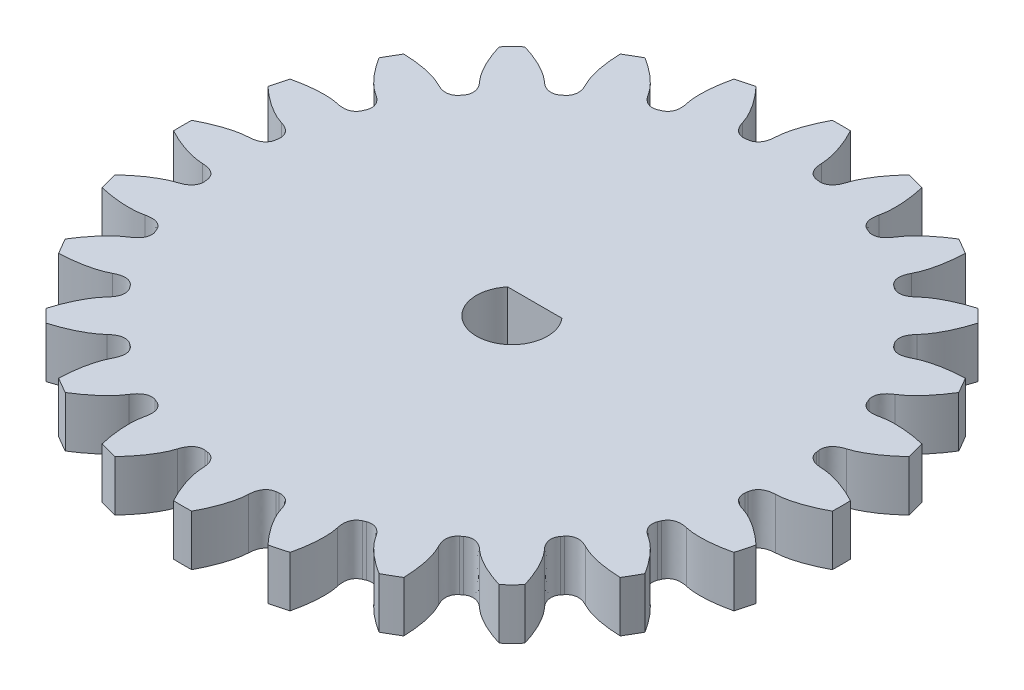
SolidWorks part; units mm, degrees
ref_plane "Спереди" through (0, 0, 0) normal (0, 0, 1) x (1, 0, 0)
ref_plane "Сверху" through (0, 0, 0) normal (0, 1, 0) x (1, 0, 0)
ref_plane "Справа" through (0, 0, 0) normal (1, 0, 0) x (0, 0, -1)
sketch "Эскиз1" plane through (0, 0, 0) normal (0, 1, 0) x (1, 0, 0)
  line L0 (-1.0724, 0.9) -> (1.0724, 0.9)
  arc A3 (-1.0724, 0.9) -> (1.0724, 0.9) centre (0, 0) ccw
  point P1 (0, -1.4)
  line B0 (-14.3, 0) -> (14.3, 0) construction
  line B1 (0, -14.3) -> (0, 14.3) construction
  arc B2 (0.3577, 12.9951) -> (-0.3577, 12.9951) centre (0, 0) ccw
  arc B3 (-1.346, 10.6654) -> (-1.4603, 10.6504) centre (0, 0) ccw
  arc B4 (-3.0178, 12.6449) -> (-3.7089, 12.4597) centre (0, 0) ccw
  arc B5 (-4.0605, 9.9536) -> (-4.1671, 9.9095) centre (0, 0) ccw
  arc B6 (-6.1877, 11.4329) -> (-6.8073, 11.0752) centre (0, 0) ccw
  arc B7 (-6.4984, 8.5635) -> (-6.5898, 8.4933) centre (0, 0) ccw
  arc B8 (-8.936, 9.4419) -> (-9.4419, 8.936) centre (0, 0) ccw
  arc B9 (-8.4933, 6.5898) -> (-8.5635, 6.4984) centre (0, 0) ccw
  arc B10 (-11.0752, 6.8073) -> (-11.4329, 6.1877) centre (0, 0) ccw
  arc B11 (-9.9095, 4.1671) -> (-9.9536, 4.0605) centre (0, 0) ccw
  arc B12 (-12.4597, 3.7089) -> (-12.6449, 3.0178) centre (0, 0) ccw
  arc B13 (-10.6504, 1.4603) -> (-10.6654, 1.346) centre (0, 0) ccw
  arc B14 (-12.9951, 0.3577) -> (-12.9951, -0.3577) centre (0, 0) ccw
  arc B15 (-10.6654, -1.346) -> (-10.6504, -1.4603) centre (0, 0) ccw
  arc B16 (-12.6449, -3.0178) -> (-12.4597, -3.7089) centre (0, 0) ccw
  arc B17 (-9.9536, -4.0605) -> (-9.9095, -4.1671) centre (0, 0) ccw
  arc B18 (-11.4329, -6.1877) -> (-11.0752, -6.8073) centre (0, 0) ccw
  arc B19 (-8.5635, -6.4984) -> (-8.4933, -6.5898) centre (0, 0) ccw
  arc B20 (-9.4419, -8.936) -> (-8.936, -9.4419) centre (0, 0) ccw
  arc B21 (-6.5898, -8.4933) -> (-6.4984, -8.5635) centre (0, 0) ccw
  arc B22 (-6.8073, -11.0752) -> (-6.1877, -11.4329) centre (0, 0) ccw
  arc B23 (-4.1671, -9.9095) -> (-4.0605, -9.9536) centre (0, 0) ccw
  arc B24 (-3.7089, -12.4597) -> (-3.0178, -12.6449) centre (0, 0) ccw
  arc B25 (-1.4603, -10.6504) -> (-1.346, -10.6654) centre (0, 0) ccw
  arc B26 (-0.3577, -12.9951) -> (0.3577, -12.9951) centre (0, 0) ccw
  arc B27 (1.346, -10.6654) -> (1.4603, -10.6504) centre (0, 0) ccw
  arc B28 (3.0178, -12.6449) -> (3.7089, -12.4597) centre (0, 0) ccw
  arc B29 (4.0605, -9.9536) -> (4.1671, -9.9095) centre (0, 0) ccw
  arc B30 (6.1877, -11.4329) -> (6.8073, -11.0752) centre (0, 0) ccw
  arc B31 (6.4984, -8.5635) -> (6.5898, -8.4933) centre (0, 0) ccw
  arc B32 (8.936, -9.4419) -> (9.4419, -8.936) centre (0, 0) ccw
  arc B33 (8.4933, -6.5898) -> (8.5635, -6.4984) centre (0, 0) ccw
  arc B34 (11.0752, -6.8073) -> (11.4329, -6.1877) centre (0, 0) ccw
  arc B35 (9.9095, -4.1671) -> (9.9536, -4.0605) centre (0, 0) ccw
  arc B36 (12.4597, -3.7089) -> (12.6449, -3.0178) centre (0, 0) ccw
  arc B37 (10.6504, -1.4603) -> (10.6654, -1.346) centre (0, 0) ccw
  arc B38 (12.9951, -0.3577) -> (12.9951, 0.3577) centre (0, 0) ccw
  arc B39 (10.6654, 1.346) -> (10.6504, 1.4603) centre (0, 0) ccw
  arc B40 (12.6449, 3.0178) -> (12.4597, 3.7089) centre (0, 0) ccw
  arc B41 (9.9536, 4.0605) -> (9.9095, 4.1671) centre (0, 0) ccw
  arc B42 (11.4329, 6.1877) -> (11.0752, 6.8073) centre (0, 0) ccw
  arc B43 (8.5635, 6.4984) -> (8.4933, 6.5898) centre (0, 0) ccw
  arc B44 (9.4419, 8.936) -> (8.936, 9.4419) centre (0, 0) ccw
  arc B45 (6.5898, 8.4933) -> (6.4984, 8.5635) centre (0, 0) ccw
  arc B46 (6.8073, 11.0752) -> (6.1877, 11.4329) centre (0, 0) ccw
  arc B47 (4.1671, 9.9095) -> (4.0605, 9.9536) centre (0, 0) ccw
  arc B48 (3.7089, 12.4597) -> (3.0178, 12.6449) centre (0, 0) ccw
  arc B49 (1.4603, 10.6504) -> (1.346, 10.6654) centre (0, 0) ccw
  circle B50 centre (0, 0) radius 12 construction
  spline B51 degree 3 poles (0.9058, 11.3017) (0.9058, 11.2304) (0.9138, 11.1608) (0.9299, 11.0929) (0.9396, 11.0522) (0.9513, 11.0113) (0.9676, 10.9727) (0.9799, 10.9437) (0.994, 10.915) (1.0107, 10.8883) (1.0248, 10.8656) (1.0406, 10.8436) (1.058, 10.8234) (1.0738, 10.805) (1.091, 10.7875) (1.1093, 10.7717) (1.1266, 10.7569) (1.1451, 10.7431) (1.1643, 10.7309) (1.1829, 10.7192) (1.2025, 10.7087) (1.2225, 10.6998) (1.2421, 10.6911) (1.2626, 10.6838) (1.2833, 10.678) (1.3038, 10.6723) (1.3247, 10.6681) (1.346, 10.6654) knots 0 0 0 0 1 1 1 2 2 2 3 3 3 4 4 4 5 5 5 6 6 6 7 7 7 8 8 8 9 9 9 9
  spline B52 degree 3 poles (-0.9058, 11.3017) (-0.9058, 11.2304) (-0.9138, 11.1608) (-0.9299, 11.0929) (-0.9396, 11.0522) (-0.9513, 11.0113) (-0.9676, 10.9727) (-0.9799, 10.9437) (-0.994, 10.915) (-1.0107, 10.8883) (-1.0248, 10.8656) (-1.0406, 10.8436) (-1.058, 10.8234) (-1.0738, 10.805) (-1.091, 10.7875) (-1.1093, 10.7717) (-1.1266, 10.7569) (-1.1451, 10.7431) (-1.1643, 10.7309) (-1.1829, 10.7192) (-1.2025, 10.7087) (-1.2225, 10.6998) (-1.2421, 10.6911) (-1.2626, 10.6838) (-1.2833, 10.678) (-1.3038, 10.6723) (-1.3247, 10.6681) (-1.346, 10.6654) knots 0 0 0 0 1 1 1 2 2 2 3 3 3 4 4 4 5 5 5 6 6 6 7 7 7 8 8 8 9 9 9 9
  spline B53 degree 3 poles (0.9058, 11.3017) (0.9032, 11.3642) (0.898, 11.4263) (0.8903, 11.4882) (0.8824, 11.551) (0.8712, 11.6136) (0.8589, 11.6757) (0.8463, 11.7389) (0.8314, 11.8016) (0.8153, 11.864) (0.7989, 11.9273) (0.7806, 11.9902) (0.7612, 12.0526) (0.7414, 12.116) (0.72, 12.179) (0.6975, 12.2415) (0.6746, 12.3049) (0.6503, 12.3678) (0.6249, 12.4303) (0.5991, 12.4937) (0.572, 12.5566) (0.5439, 12.6189) (0.5153, 12.6822) (0.4855, 12.745) (0.4547, 12.8073) (0.4235, 12.8704) (0.3912, 12.933) (0.3577, 12.9951) knots 0 0 0 0 1 1 1 2 2 2 3 3 3 4 4 4 5 5 5 6 6 6 7 7 7 8 8 8 9 9 9 9
  spline B54 degree 3 poles (-0.9058, 11.3017) (-0.9032, 11.3642) (-0.898, 11.4263) (-0.8903, 11.4882) (-0.8824, 11.551) (-0.8712, 11.6136) (-0.8589, 11.6757) (-0.8463, 11.7389) (-0.8314, 11.8016) (-0.8153, 11.864) (-0.7989, 11.9273) (-0.7806, 11.9902) (-0.7612, 12.0526) (-0.7414, 12.116) (-0.72, 12.179) (-0.6975, 12.2415) (-0.6746, 12.3049) (-0.6503, 12.3678) (-0.6249, 12.4303) (-0.5991, 12.4937) (-0.572, 12.5566) (-0.5439, 12.6189) (-0.5153, 12.6822) (-0.4855, 12.745) (-0.4547, 12.8073) (-0.4235, 12.8704) (-0.3912, 12.933) (-0.3577, 12.9951) knots 0 0 0 0 1 1 1 2 2 2 3 3 3 4 4 4 5 5 5 6 6 6 7 7 7 8 8 8 9 9 9 9
  spline B55 degree 3 poles (-2.0502, 11.151) (-2.0317, 11.0822) (-2.0059, 11.017) (-1.9728, 10.9556) (-1.9529, 10.9188) (-1.931, 10.8823) (-1.9053, 10.8493) (-1.886, 10.8244) (-1.8649, 10.8004) (-1.8419, 10.7789) (-1.8224, 10.7606) (-1.8014, 10.7435) (-1.7793, 10.7284) (-1.7594, 10.7148) (-1.7382, 10.7023) (-1.7164, 10.6918) (-1.6959, 10.6819) (-1.6745, 10.6734) (-1.6527, 10.6666) (-1.6318, 10.6601) (-1.6101, 10.655) (-1.5885, 10.6516) (-1.5672, 10.6483) (-1.5456, 10.6465) (-1.5241, 10.6463) (-1.5028, 10.6461) (-1.4816, 10.6475) (-1.4603, 10.6504) knots 0 0 0 0 1 1 1 2 2 2 3 3 3 4 4 4 5 5 5 6 6 6 7 7 7 8 8 8 9 9 9 9
  spline B56 degree 3 poles (-3.8, 10.6822) (-3.7815, 10.6133) (-3.7713, 10.544) (-3.7693, 10.4743) (-3.7681, 10.4325) (-3.7688, 10.3898) (-3.7746, 10.3484) (-3.7789, 10.3172) (-3.7852, 10.2858) (-3.7943, 10.2557) (-3.8021, 10.2302) (-3.8117, 10.2048) (-3.8232, 10.1807) (-3.8337, 10.1589) (-3.8458, 10.1376) (-3.8595, 10.1176) (-3.8723, 10.0988) (-3.8866, 10.0806) (-3.902, 10.0639) (-3.9169, 10.0478) (-3.9331, 10.0326) (-3.9502, 10.0188) (-3.9669, 10.0053) (-3.9848, 9.9929) (-4.0032, 9.982) (-4.0216, 9.9712) (-4.0406, 9.9618) (-4.0605, 9.9536) knots 0 0 0 0 1 1 1 2 2 2 3 3 3 4 4 4 5 5 5 6 6 6 7 7 7 8 8 8 9 9 9 9
  spline B57 degree 3 poles (-2.0502, 11.151) (-2.0689, 11.2107) (-2.09, 11.2694) (-2.1134, 11.3271) (-2.1373, 11.3858) (-2.1643, 11.4434) (-2.1923, 11.5002) (-2.2208, 11.5579) (-2.2514, 11.6147) (-2.2831, 11.6707) (-2.3153, 11.7276) (-2.3493, 11.7837) (-2.3842, 11.8389) (-2.4197, 11.8951) (-2.4567, 11.9503) (-2.4946, 12.0049) (-2.5331, 12.0602) (-2.5729, 12.1147) (-2.6136, 12.1685) (-2.6549, 12.223) (-2.6974, 12.2768) (-2.7407, 12.3297) (-2.7847, 12.3835) (-2.8297, 12.4364) (-2.8755, 12.4885) (-2.9221, 12.5415) (-2.9695, 12.5936) (-3.0178, 12.6449) knots 0 0 0 0 1 1 1 2 2 2 3 3 3 4 4 4 5 5 5 6 6 6 7 7 7 8 8 8 9 9 9 9
  spline B58 degree 3 poles (-3.8, 10.6822) (-3.8136, 10.7432) (-3.8247, 10.8046) (-3.8333, 10.8663) (-3.842, 10.929) (-3.8474, 10.9924) (-3.8515, 11.0556) (-3.8557, 11.1198) (-3.8576, 11.1843) (-3.8581, 11.2487) (-3.8587, 11.3141) (-3.8573, 11.3796) (-3.8547, 11.4449) (-3.852, 11.5113) (-3.8476, 11.5776) (-3.8421, 11.6438) (-3.8364, 11.711) (-3.8292, 11.7781) (-3.8208, 11.845) (-3.8123, 11.9129) (-3.8024, 11.9807) (-3.7914, 12.0482) (-3.7802, 12.1167) (-3.7676, 12.1851) (-3.754, 12.2532) (-3.7402, 12.3223) (-3.7251, 12.3911) (-3.7089, 12.4597) knots 0 0 0 0 1 1 1 2 2 2 3 3 3 4 4 4 5 5 5 6 6 6 7 7 7 8 8 8 9 9 9 9
  spline B59 degree 3 poles (-4.8664, 10.2404) (-4.8308, 10.1787) (-4.789, 10.1225) (-4.7411, 10.0717) (-4.7124, 10.0413) (-4.6817, 10.0117) (-4.6484, 9.9865) (-4.6233, 9.9675) (-4.5967, 9.9497) (-4.5689, 9.9349) (-4.5453, 9.9223) (-4.5206, 9.9111) (-4.4954, 9.9023) (-4.4726, 9.8943) (-4.4489, 9.8878) (-4.4252, 9.8833) (-4.4028, 9.879) (-4.3799, 9.8763) (-4.3571, 9.8754) (-4.3352, 9.8745) (-4.313, 9.8752) (-4.2912, 9.8776) (-4.2698, 9.8798) (-4.2484, 9.8837) (-4.2276, 9.8891) (-4.2071, 9.8944) (-4.1869, 9.9012) (-4.1671, 9.9095) knots 0 0 0 0 1 1 1 2 2 2 3 3 3 4 4 4 5 5 5 6 6 6 7 7 7 8 8 8 9 9 9 9
  spline B60 degree 3 poles (-6.4353, 9.3347) (-6.3996, 9.2729) (-6.3718, 9.2086) (-6.3518, 9.1418) (-6.3398, 9.1017) (-6.3295, 9.0604) (-6.3243, 9.0188) (-6.3204, 8.9876) (-6.3184, 8.9557) (-6.3194, 8.9242) (-6.3203, 8.8975) (-6.323, 8.8706) (-6.3279, 8.8443) (-6.3324, 8.8205) (-6.3386, 8.7968) (-6.3466, 8.7739) (-6.3541, 8.7524) (-6.3632, 8.7312) (-6.3738, 8.7111) (-6.384, 8.6917) (-6.3957, 8.6728) (-6.4086, 8.655) (-6.4213, 8.6377) (-6.4353, 8.6211) (-6.4504, 8.6058) (-6.4653, 8.5906) (-6.4813, 8.5765) (-6.4984, 8.5635) knots 0 0 0 0 1 1 1 2 2 2 3 3 3 4 4 4 5 5 5 6 6 6 7 7 7 8 8 8 9 9 9 9
  spline B61 degree 3 poles (-4.8664, 10.2404) (-4.8999, 10.2932) (-4.9355, 10.3445) (-4.9731, 10.3942) (-5.0113, 10.4447) (-5.0523, 10.4933) (-5.0941, 10.5409) (-5.1365, 10.5893) (-5.1808, 10.6362) (-5.2259, 10.6822) (-5.2718, 10.7288) (-5.319, 10.7741) (-5.3671, 10.8185) (-5.4159, 10.8635) (-5.4659, 10.9073) (-5.5167, 10.9502) (-5.5682, 10.9937) (-5.6207, 11.036) (-5.674, 11.0774) (-5.728, 11.1194) (-5.7829, 11.1603) (-5.8385, 11.2003) (-5.8949, 11.2408) (-5.9521, 11.2803) (-6.0098, 11.3188) (-6.0685, 11.3578) (-6.1278, 11.3959) (-6.1877, 11.4329) knots 0 0 0 0 1 1 1 2 2 2 3 3 3 4 4 4 5 5 5 6 6 6 7 7 7 8 8 8 9 9 9 9
  spline B62 degree 3 poles (-6.4353, 9.3347) (-6.4642, 9.3901) (-6.4908, 9.4465) (-6.5151, 9.5039) (-6.5397, 9.5623) (-6.5613, 9.622) (-6.5817, 9.6821) (-6.6024, 9.743) (-6.6209, 9.8048) (-6.638, 9.8669) (-6.6555, 9.9299) (-6.6711, 9.9935) (-6.6855, 10.0573) (-6.7001, 10.1221) (-6.713, 10.1873) (-6.7248, 10.2527) (-6.7367, 10.319) (-6.7471, 10.3857) (-6.7563, 10.4525) (-6.7657, 10.5203) (-6.7737, 10.5883) (-6.7805, 10.6564) (-6.7874, 10.7255) (-6.793, 10.7948) (-6.7974, 10.8641) (-6.8019, 10.9344) (-6.8053, 11.0047) (-6.8073, 11.0752) knots 0 0 0 0 1 1 1 2 2 2 3 3 3 4 4 4 5 5 5 6 6 6 7 7 7 8 8 8 9 9 9 9
  spline B63 degree 3 poles (-7.351, 8.632) (-7.3006, 8.5816) (-7.2457, 8.5381) (-7.1863, 8.5015) (-7.1507, 8.4795) (-7.1134, 8.4588) (-7.0747, 8.4431) (-7.0455, 8.4312) (-7.0152, 8.421) (-6.9845, 8.4138) (-6.9585, 8.4078) (-6.9318, 8.4034) (-6.9052, 8.4014) (-6.881, 8.3996) (-6.8565, 8.3994) (-6.8324, 8.4012) (-6.8097, 8.4029) (-6.7868, 8.4062) (-6.7646, 8.4112) (-6.7432, 8.416) (-6.7219, 8.4224) (-6.7015, 8.4304) (-6.6814, 8.4381) (-6.6618, 8.4474) (-6.6431, 8.4579) (-6.6246, 8.4684) (-6.6068, 8.4802) (-6.5898, 8.4933) knots 0 0 0 0 1 1 1 2 2 2 3 3 3 4 4 4 5 5 5 6 6 6 7 7 7 8 8 8 9 9 9 9
  spline B64 degree 3 poles (-8.632, 7.351) (-8.5816, 7.3006) (-8.5381, 7.2457) (-8.5015, 7.1863) (-8.4795, 7.1507) (-8.4588, 7.1134) (-8.4431, 7.0747) (-8.4312, 7.0455) (-8.421, 7.0152) (-8.4138, 6.9845) (-8.4078, 6.9585) (-8.4034, 6.9318) (-8.4014, 6.9052) (-8.3996, 6.881) (-8.3994, 6.8565) (-8.4012, 6.8324) (-8.4029, 6.8097) (-8.4062, 6.7868) (-8.4112, 6.7646) (-8.416, 6.7432) (-8.4224, 6.7219) (-8.4304, 6.7015) (-8.4381, 6.6814) (-8.4474, 6.6618) (-8.4579, 6.6431) (-8.4684, 6.6246) (-8.4802, 6.6068) (-8.4933, 6.5898) knots 0 0 0 0 1 1 1 2 2 2 3 3 3 4 4 4 5 5 5 6 6 6 7 7 7 8 8 8 9 9 9 9
  spline B65 degree 3 poles (-7.351, 8.632) (-7.3971, 8.6743) (-7.4447, 8.7146) (-7.4938, 8.7529) (-7.5438, 8.7918) (-7.596, 8.8281) (-7.6487, 8.8633) (-7.7022, 8.8991) (-7.7571, 8.9329) (-7.8126, 8.9656) (-7.869, 8.9988) (-7.9263, 9.0303) (-7.9843, 9.0607) (-8.0431, 9.0916) (-8.1027, 9.121) (-8.1628, 9.1492) (-8.2238, 9.1779) (-8.2855, 9.2052) (-8.3477, 9.2314) (-8.4107, 9.258) (-8.4744, 9.2833) (-8.5384, 9.3075) (-8.6033, 9.3321) (-8.6688, 9.3554) (-8.7346, 9.3776) (-8.8013, 9.4002) (-8.8684, 9.4216) (-8.936, 9.4419) knots 0 0 0 0 1 1 1 2 2 2 3 3 3 4 4 4 5 5 5 6 6 6 7 7 7 8 8 8 9 9 9 9
  spline B66 degree 3 poles (-8.632, 7.351) (-8.6743, 7.3971) (-8.7146, 7.4447) (-8.7529, 7.4938) (-8.7918, 7.5438) (-8.8281, 7.596) (-8.8633, 7.6487) (-8.8991, 7.7022) (-8.9329, 7.7571) (-8.9656, 7.8126) (-8.9988, 7.869) (-9.0303, 7.9263) (-9.0607, 7.9843) (-9.0916, 8.0431) (-9.121, 8.1027) (-9.1492, 8.1628) (-9.1779, 8.2238) (-9.2052, 8.2855) (-9.2314, 8.3477) (-9.258, 8.4107) (-9.2833, 8.4744) (-9.3075, 8.5384) (-9.3321, 8.6033) (-9.3554, 8.6688) (-9.3776, 8.7346) (-9.4002, 8.8013) (-9.4216, 8.8684) (-9.4419, 8.936) knots 0 0 0 0 1 1 1 2 2 2 3 3 3 4 4 4 5 5 5 6 6 6 7 7 7 8 8 8 9 9 9 9
  spline B67 degree 3 poles (-9.3347, 6.4353) (-9.2729, 6.3996) (-9.2086, 6.3718) (-9.1418, 6.3518) (-9.1017, 6.3398) (-9.0604, 6.3295) (-9.0188, 6.3243) (-8.9876, 6.3204) (-8.9557, 6.3184) (-8.9242, 6.3194) (-8.8975, 6.3203) (-8.8706, 6.323) (-8.8443, 6.3279) (-8.8205, 6.3324) (-8.7968, 6.3386) (-8.7739, 6.3466) (-8.7524, 6.3541) (-8.7312, 6.3632) (-8.7111, 6.3738) (-8.6917, 6.384) (-8.6728, 6.3957) (-8.655, 6.4086) (-8.6377, 6.4213) (-8.6211, 6.4353) (-8.6058, 6.4504) (-8.5906, 6.4653) (-8.5765, 6.4813) (-8.5635, 6.4984) knots 0 0 0 0 1 1 1 2 2 2 3 3 3 4 4 4 5 5 5 6 6 6 7 7 7 8 8 8 9 9 9 9
  spline B68 degree 3 poles (-10.2404, 4.8664) (-10.1787, 4.8308) (-10.1225, 4.789) (-10.0717, 4.7411) (-10.0413, 4.7124) (-10.0117, 4.6817) (-9.9865, 4.6484) (-9.9675, 4.6233) (-9.9497, 4.5967) (-9.9349, 4.5689) (-9.9223, 4.5453) (-9.9111, 4.5206) (-9.9023, 4.4954) (-9.8943, 4.4726) (-9.8878, 4.4489) (-9.8833, 4.4252) (-9.879, 4.4028) (-9.8763, 4.3799) (-9.8754, 4.3571) (-9.8745, 4.3352) (-9.8752, 4.313) (-9.8776, 4.2912) (-9.8798, 4.2698) (-9.8837, 4.2484) (-9.8891, 4.2276) (-9.8944, 4.2071) (-9.9012, 4.1869) (-9.9095, 4.1671) knots 0 0 0 0 1 1 1 2 2 2 3 3 3 4 4 4 5 5 5 6 6 6 7 7 7 8 8 8 9 9 9 9
  spline B69 degree 3 poles (-9.3347, 6.4353) (-9.3901, 6.4642) (-9.4465, 6.4908) (-9.5039, 6.5151) (-9.5623, 6.5397) (-9.622, 6.5613) (-9.6821, 6.5817) (-9.743, 6.6024) (-9.8048, 6.6209) (-9.8669, 6.638) (-9.9299, 6.6555) (-9.9935, 6.6711) (-10.0573, 6.6855) (-10.1221, 6.7001) (-10.1873, 6.713) (-10.2527, 6.7248) (-10.319, 6.7367) (-10.3857, 6.7471) (-10.4525, 6.7563) (-10.5203, 6.7657) (-10.5883, 6.7737) (-10.6564, 6.7805) (-10.7255, 6.7874) (-10.7948, 6.793) (-10.8641, 6.7974) (-10.9344, 6.8019) (-11.0047, 6.8053) (-11.0752, 6.8073) knots 0 0 0 0 1 1 1 2 2 2 3 3 3 4 4 4 5 5 5 6 6 6 7 7 7 8 8 8 9 9 9 9
  spline B70 degree 3 poles (-10.2404, 4.8664) (-10.2932, 4.8999) (-10.3445, 4.9355) (-10.3942, 4.9731) (-10.4447, 5.0113) (-10.4933, 5.0523) (-10.5409, 5.0941) (-10.5893, 5.1365) (-10.6362, 5.1808) (-10.6822, 5.2259) (-10.7288, 5.2718) (-10.7741, 5.319) (-10.8185, 5.3671) (-10.8635, 5.4159) (-10.9073, 5.4659) (-10.9502, 5.5167) (-10.9937, 5.5682) (-11.036, 5.6207) (-11.0774, 5.674) (-11.1194, 5.728) (-11.1603, 5.7829) (-11.2003, 5.8385) (-11.2408, 5.8949) (-11.2803, 5.9521) (-11.3188, 6.0098) (-11.3578, 6.0685) (-11.3959, 6.1278) (-11.4329, 6.1877) knots 0 0 0 0 1 1 1 2 2 2 3 3 3 4 4 4 5 5 5 6 6 6 7 7 7 8 8 8 9 9 9 9
  spline B71 degree 3 poles (-10.6822, 3.8) (-10.6133, 3.7815) (-10.544, 3.7713) (-10.4743, 3.7693) (-10.4325, 3.7681) (-10.3898, 3.7688) (-10.3484, 3.7746) (-10.3172, 3.7789) (-10.2858, 3.7852) (-10.2557, 3.7943) (-10.2302, 3.8021) (-10.2048, 3.8117) (-10.1807, 3.8232) (-10.1589, 3.8337) (-10.1376, 3.8458) (-10.1176, 3.8595) (-10.0988, 3.8723) (-10.0806, 3.8866) (-10.0639, 3.902) (-10.0478, 3.9169) (-10.0326, 3.9331) (-10.0188, 3.9502) (-10.0053, 3.9669) (-9.9929, 3.9848) (-9.982, 4.0032) (-9.9712, 4.0216) (-9.9618, 4.0406) (-9.9536, 4.0605) knots 0 0 0 0 1 1 1 2 2 2 3 3 3 4 4 4 5 5 5 6 6 6 7 7 7 8 8 8 9 9 9 9
  spline B72 degree 3 poles (-11.151, 2.0502) (-11.0822, 2.0317) (-11.017, 2.0059) (-10.9556, 1.9728) (-10.9188, 1.9529) (-10.8823, 1.931) (-10.8493, 1.9053) (-10.8244, 1.886) (-10.8004, 1.8649) (-10.7789, 1.8419) (-10.7606, 1.8224) (-10.7435, 1.8014) (-10.7284, 1.7793) (-10.7148, 1.7594) (-10.7023, 1.7382) (-10.6918, 1.7164) (-10.6819, 1.6959) (-10.6734, 1.6745) (-10.6666, 1.6527) (-10.6601, 1.6318) (-10.655, 1.6101) (-10.6516, 1.5885) (-10.6483, 1.5672) (-10.6465, 1.5456) (-10.6463, 1.5241) (-10.6461, 1.5028) (-10.6475, 1.4816) (-10.6504, 1.4603) knots 0 0 0 0 1 1 1 2 2 2 3 3 3 4 4 4 5 5 5 6 6 6 7 7 7 8 8 8 9 9 9 9
  spline B73 degree 3 poles (-10.6822, 3.8) (-10.7432, 3.8136) (-10.8046, 3.8247) (-10.8663, 3.8333) (-10.929, 3.842) (-10.9924, 3.8474) (-11.0556, 3.8515) (-11.1198, 3.8557) (-11.1843, 3.8576) (-11.2487, 3.8581) (-11.3141, 3.8587) (-11.3796, 3.8573) (-11.4449, 3.8547) (-11.5113, 3.852) (-11.5776, 3.8476) (-11.6438, 3.8421) (-11.711, 3.8364) (-11.7781, 3.8292) (-11.845, 3.8208) (-11.9129, 3.8123) (-11.9807, 3.8024) (-12.0482, 3.7914) (-12.1167, 3.7802) (-12.1851, 3.7676) (-12.2532, 3.754) (-12.3223, 3.7402) (-12.3911, 3.7251) (-12.4597, 3.7089) knots 0 0 0 0 1 1 1 2 2 2 3 3 3 4 4 4 5 5 5 6 6 6 7 7 7 8 8 8 9 9 9 9
  spline B74 degree 3 poles (-11.151, 2.0502) (-11.2107, 2.0689) (-11.2694, 2.09) (-11.3271, 2.1134) (-11.3858, 2.1373) (-11.4434, 2.1643) (-11.5002, 2.1923) (-11.5579, 2.2208) (-11.6147, 2.2514) (-11.6707, 2.2831) (-11.7276, 2.3153) (-11.7837, 2.3493) (-11.8389, 2.3842) (-11.8951, 2.4197) (-11.9503, 2.4567) (-12.0049, 2.4946) (-12.0602, 2.5331) (-12.1147, 2.5729) (-12.1685, 2.6136) (-12.223, 2.6549) (-12.2768, 2.6974) (-12.3297, 2.7407) (-12.3835, 2.7847) (-12.4364, 2.8297) (-12.4885, 2.8755) (-12.5415, 2.9221) (-12.5936, 2.9695) (-12.6449, 3.0178) knots 0 0 0 0 1 1 1 2 2 2 3 3 3 4 4 4 5 5 5 6 6 6 7 7 7 8 8 8 9 9 9 9
  spline B75 degree 3 poles (-11.3017, 0.9058) (-11.2304, 0.9058) (-11.1608, 0.9138) (-11.0929, 0.9299) (-11.0522, 0.9396) (-11.0113, 0.9513) (-10.9727, 0.9676) (-10.9437, 0.9799) (-10.915, 0.994) (-10.8883, 1.0107) (-10.8656, 1.0248) (-10.8436, 1.0406) (-10.8234, 1.058) (-10.805, 1.0738) (-10.7875, 1.091) (-10.7717, 1.1093) (-10.7569, 1.1266) (-10.7431, 1.1451) (-10.7309, 1.1643) (-10.7192, 1.1829) (-10.7087, 1.2025) (-10.6998, 1.2225) (-10.6911, 1.2421) (-10.6838, 1.2626) (-10.678, 1.2833) (-10.6723, 1.3038) (-10.6681, 1.3247) (-10.6654, 1.346) knots 0 0 0 0 1 1 1 2 2 2 3 3 3 4 4 4 5 5 5 6 6 6 7 7 7 8 8 8 9 9 9 9
  spline B76 degree 3 poles (-11.3017, -0.9058) (-11.2304, -0.9058) (-11.1608, -0.9138) (-11.0929, -0.9299) (-11.0522, -0.9396) (-11.0113, -0.9513) (-10.9727, -0.9676) (-10.9437, -0.9799) (-10.915, -0.994) (-10.8883, -1.0107) (-10.8656, -1.0248) (-10.8436, -1.0406) (-10.8234, -1.058) (-10.805, -1.0738) (-10.7875, -1.091) (-10.7717, -1.1093) (-10.7569, -1.1266) (-10.7431, -1.1451) (-10.7309, -1.1643) (-10.7192, -1.1829) (-10.7087, -1.2025) (-10.6998, -1.2225) (-10.6911, -1.2421) (-10.6838, -1.2626) (-10.678, -1.2833) (-10.6723, -1.3038) (-10.6681, -1.3247) (-10.6654, -1.346) knots 0 0 0 0 1 1 1 2 2 2 3 3 3 4 4 4 5 5 5 6 6 6 7 7 7 8 8 8 9 9 9 9
  spline B77 degree 3 poles (-11.3017, 0.9058) (-11.3642, 0.9032) (-11.4263, 0.898) (-11.4882, 0.8903) (-11.551, 0.8824) (-11.6136, 0.8712) (-11.6757, 0.8589) (-11.7389, 0.8463) (-11.8016, 0.8314) (-11.864, 0.8153) (-11.9273, 0.7989) (-11.9902, 0.7806) (-12.0526, 0.7612) (-12.116, 0.7414) (-12.179, 0.72) (-12.2415, 0.6975) (-12.3049, 0.6746) (-12.3678, 0.6503) (-12.4303, 0.6249) (-12.4937, 0.5991) (-12.5566, 0.572) (-12.6189, 0.5439) (-12.6822, 0.5153) (-12.745, 0.4855) (-12.8073, 0.4547) (-12.8704, 0.4235) (-12.933, 0.3912) (-12.9951, 0.3577) knots 0 0 0 0 1 1 1 2 2 2 3 3 3 4 4 4 5 5 5 6 6 6 7 7 7 8 8 8 9 9 9 9
  spline B78 degree 3 poles (-11.3017, -0.9058) (-11.3642, -0.9032) (-11.4263, -0.898) (-11.4882, -0.8903) (-11.551, -0.8824) (-11.6136, -0.8712) (-11.6757, -0.8589) (-11.7389, -0.8463) (-11.8016, -0.8314) (-11.864, -0.8153) (-11.9273, -0.7989) (-11.9902, -0.7806) (-12.0526, -0.7612) (-12.116, -0.7414) (-12.179, -0.72) (-12.2415, -0.6975) (-12.3049, -0.6746) (-12.3678, -0.6503) (-12.4303, -0.6249) (-12.4937, -0.5991) (-12.5566, -0.572) (-12.6189, -0.5439) (-12.6822, -0.5153) (-12.745, -0.4855) (-12.8073, -0.4547) (-12.8704, -0.4235) (-12.933, -0.3912) (-12.9951, -0.3577) knots 0 0 0 0 1 1 1 2 2 2 3 3 3 4 4 4 5 5 5 6 6 6 7 7 7 8 8 8 9 9 9 9
  spline B79 degree 3 poles (-11.151, -2.0502) (-11.0822, -2.0317) (-11.017, -2.0059) (-10.9556, -1.9728) (-10.9188, -1.9529) (-10.8823, -1.931) (-10.8493, -1.9053) (-10.8244, -1.886) (-10.8004, -1.8649) (-10.7789, -1.8419) (-10.7606, -1.8224) (-10.7435, -1.8014) (-10.7284, -1.7793) (-10.7148, -1.7594) (-10.7023, -1.7382) (-10.6918, -1.7164) (-10.6819, -1.6959) (-10.6734, -1.6745) (-10.6666, -1.6527) (-10.6601, -1.6318) (-10.655, -1.6101) (-10.6516, -1.5885) (-10.6483, -1.5672) (-10.6465, -1.5456) (-10.6463, -1.5241) (-10.6461, -1.5028) (-10.6475, -1.4816) (-10.6504, -1.4603) knots 0 0 0 0 1 1 1 2 2 2 3 3 3 4 4 4 5 5 5 6 6 6 7 7 7 8 8 8 9 9 9 9
  spline B80 degree 3 poles (-10.6822, -3.8) (-10.6133, -3.7815) (-10.544, -3.7713) (-10.4743, -3.7693) (-10.4325, -3.7681) (-10.3898, -3.7688) (-10.3484, -3.7746) (-10.3172, -3.7789) (-10.2858, -3.7852) (-10.2557, -3.7943) (-10.2302, -3.8021) (-10.2048, -3.8117) (-10.1807, -3.8232) (-10.1589, -3.8337) (-10.1376, -3.8458) (-10.1176, -3.8595) (-10.0988, -3.8723) (-10.0806, -3.8866) (-10.0639, -3.902) (-10.0478, -3.9169) (-10.0326, -3.9331) (-10.0188, -3.9502) (-10.0053, -3.9669) (-9.9929, -3.9848) (-9.982, -4.0032) (-9.9712, -4.0216) (-9.9618, -4.0406) (-9.9536, -4.0605) knots 0 0 0 0 1 1 1 2 2 2 3 3 3 4 4 4 5 5 5 6 6 6 7 7 7 8 8 8 9 9 9 9
  spline B81 degree 3 poles (-11.151, -2.0502) (-11.2107, -2.0689) (-11.2694, -2.09) (-11.3271, -2.1134) (-11.3858, -2.1373) (-11.4434, -2.1643) (-11.5002, -2.1923) (-11.5579, -2.2208) (-11.6147, -2.2514) (-11.6707, -2.2831) (-11.7276, -2.3153) (-11.7837, -2.3493) (-11.8389, -2.3842) (-11.8951, -2.4197) (-11.9503, -2.4567) (-12.0049, -2.4946) (-12.0602, -2.5331) (-12.1147, -2.5729) (-12.1685, -2.6136) (-12.223, -2.6549) (-12.2768, -2.6974) (-12.3297, -2.7407) (-12.3835, -2.7847) (-12.4364, -2.8297) (-12.4885, -2.8755) (-12.5415, -2.9221) (-12.5936, -2.9695) (-12.6449, -3.0178) knots 0 0 0 0 1 1 1 2 2 2 3 3 3 4 4 4 5 5 5 6 6 6 7 7 7 8 8 8 9 9 9 9
  spline B82 degree 3 poles (-10.6822, -3.8) (-10.7432, -3.8136) (-10.8046, -3.8247) (-10.8663, -3.8333) (-10.929, -3.842) (-10.9924, -3.8474) (-11.0556, -3.8515) (-11.1198, -3.8557) (-11.1843, -3.8576) (-11.2487, -3.8581) (-11.3141, -3.8587) (-11.3796, -3.8573) (-11.4449, -3.8547) (-11.5113, -3.852) (-11.5776, -3.8476) (-11.6438, -3.8421) (-11.711, -3.8364) (-11.7781, -3.8292) (-11.845, -3.8208) (-11.9129, -3.8123) (-11.9807, -3.8024) (-12.0482, -3.7914) (-12.1167, -3.7802) (-12.1851, -3.7676) (-12.2532, -3.754) (-12.3223, -3.7402) (-12.3911, -3.7251) (-12.4597, -3.7089) knots 0 0 0 0 1 1 1 2 2 2 3 3 3 4 4 4 5 5 5 6 6 6 7 7 7 8 8 8 9 9 9 9
  spline B83 degree 3 poles (-10.2404, -4.8664) (-10.1787, -4.8308) (-10.1225, -4.789) (-10.0717, -4.7411) (-10.0413, -4.7124) (-10.0117, -4.6817) (-9.9865, -4.6484) (-9.9675, -4.6233) (-9.9497, -4.5967) (-9.9349, -4.5689) (-9.9223, -4.5453) (-9.9111, -4.5206) (-9.9023, -4.4954) (-9.8943, -4.4726) (-9.8878, -4.4489) (-9.8833, -4.4252) (-9.879, -4.4028) (-9.8763, -4.3799) (-9.8754, -4.3571) (-9.8745, -4.3352) (-9.8752, -4.313) (-9.8776, -4.2912) (-9.8798, -4.2698) (-9.8837, -4.2484) (-9.8891, -4.2276) (-9.8944, -4.2071) (-9.9012, -4.1869) (-9.9095, -4.1671) knots 0 0 0 0 1 1 1 2 2 2 3 3 3 4 4 4 5 5 5 6 6 6 7 7 7 8 8 8 9 9 9 9
  spline B84 degree 3 poles (-9.3347, -6.4353) (-9.2729, -6.3996) (-9.2086, -6.3718) (-9.1418, -6.3518) (-9.1017, -6.3398) (-9.0604, -6.3295) (-9.0188, -6.3243) (-8.9876, -6.3204) (-8.9557, -6.3184) (-8.9242, -6.3194) (-8.8975, -6.3203) (-8.8706, -6.323) (-8.8443, -6.3279) (-8.8205, -6.3324) (-8.7968, -6.3386) (-8.7739, -6.3466) (-8.7524, -6.3541) (-8.7312, -6.3632) (-8.7111, -6.3738) (-8.6917, -6.384) (-8.6728, -6.3957) (-8.655, -6.4086) (-8.6377, -6.4213) (-8.6211, -6.4353) (-8.6058, -6.4504) (-8.5906, -6.4653) (-8.5765, -6.4813) (-8.5635, -6.4984) knots 0 0 0 0 1 1 1 2 2 2 3 3 3 4 4 4 5 5 5 6 6 6 7 7 7 8 8 8 9 9 9 9
  spline B85 degree 3 poles (-10.2404, -4.8664) (-10.2932, -4.8999) (-10.3445, -4.9355) (-10.3942, -4.9731) (-10.4447, -5.0113) (-10.4933, -5.0523) (-10.5409, -5.0941) (-10.5893, -5.1365) (-10.6362, -5.1808) (-10.6822, -5.2259) (-10.7288, -5.2718) (-10.7741, -5.319) (-10.8185, -5.3671) (-10.8635, -5.4159) (-10.9073, -5.4659) (-10.9502, -5.5167) (-10.9937, -5.5682) (-11.036, -5.6207) (-11.0774, -5.674) (-11.1194, -5.728) (-11.1603, -5.7829) (-11.2003, -5.8385) (-11.2408, -5.8949) (-11.2803, -5.9521) (-11.3188, -6.0098) (-11.3578, -6.0685) (-11.3959, -6.1278) (-11.4329, -6.1877) knots 0 0 0 0 1 1 1 2 2 2 3 3 3 4 4 4 5 5 5 6 6 6 7 7 7 8 8 8 9 9 9 9
  spline B86 degree 3 poles (-9.3347, -6.4353) (-9.3901, -6.4642) (-9.4465, -6.4908) (-9.5039, -6.5151) (-9.5623, -6.5397) (-9.622, -6.5613) (-9.6821, -6.5817) (-9.743, -6.6024) (-9.8048, -6.6209) (-9.8669, -6.638) (-9.9299, -6.6555) (-9.9935, -6.6711) (-10.0573, -6.6855) (-10.1221, -6.7001) (-10.1873, -6.713) (-10.2527, -6.7248) (-10.319, -6.7367) (-10.3857, -6.7471) (-10.4525, -6.7563) (-10.5203, -6.7657) (-10.5883, -6.7737) (-10.6564, -6.7805) (-10.7255, -6.7874) (-10.7948, -6.793) (-10.8641, -6.7974) (-10.9344, -6.8019) (-11.0047, -6.8053) (-11.0752, -6.8073) knots 0 0 0 0 1 1 1 2 2 2 3 3 3 4 4 4 5 5 5 6 6 6 7 7 7 8 8 8 9 9 9 9
  spline B87 degree 3 poles (-8.632, -7.351) (-8.5816, -7.3006) (-8.5381, -7.2457) (-8.5015, -7.1863) (-8.4795, -7.1507) (-8.4588, -7.1134) (-8.4431, -7.0747) (-8.4312, -7.0455) (-8.421, -7.0152) (-8.4138, -6.9845) (-8.4078, -6.9585) (-8.4034, -6.9318) (-8.4014, -6.9052) (-8.3996, -6.881) (-8.3994, -6.8565) (-8.4012, -6.8324) (-8.4029, -6.8097) (-8.4062, -6.7868) (-8.4112, -6.7646) (-8.416, -6.7432) (-8.4224, -6.7219) (-8.4304, -6.7015) (-8.4381, -6.6814) (-8.4474, -6.6618) (-8.4579, -6.6431) (-8.4684, -6.6246) (-8.4802, -6.6068) (-8.4933, -6.5898) knots 0 0 0 0 1 1 1 2 2 2 3 3 3 4 4 4 5 5 5 6 6 6 7 7 7 8 8 8 9 9 9 9
  spline B88 degree 3 poles (-7.351, -8.632) (-7.3006, -8.5816) (-7.2457, -8.5381) (-7.1863, -8.5015) (-7.1507, -8.4795) (-7.1134, -8.4588) (-7.0747, -8.4431) (-7.0455, -8.4312) (-7.0152, -8.421) (-6.9845, -8.4138) (-6.9585, -8.4078) (-6.9318, -8.4034) (-6.9052, -8.4014) (-6.881, -8.3996) (-6.8565, -8.3994) (-6.8324, -8.4012) (-6.8097, -8.4029) (-6.7868, -8.4062) (-6.7646, -8.4112) (-6.7432, -8.416) (-6.7219, -8.4224) (-6.7015, -8.4304) (-6.6814, -8.4381) (-6.6618, -8.4474) (-6.6431, -8.4579) (-6.6246, -8.4684) (-6.6068, -8.4802) (-6.5898, -8.4933) knots 0 0 0 0 1 1 1 2 2 2 3 3 3 4 4 4 5 5 5 6 6 6 7 7 7 8 8 8 9 9 9 9
  spline B89 degree 3 poles (-8.632, -7.351) (-8.6743, -7.3971) (-8.7146, -7.4447) (-8.7529, -7.4938) (-8.7918, -7.5438) (-8.8281, -7.596) (-8.8633, -7.6487) (-8.8991, -7.7022) (-8.9329, -7.7571) (-8.9656, -7.8126) (-8.9988, -7.869) (-9.0303, -7.9263) (-9.0607, -7.9843) (-9.0916, -8.0431) (-9.121, -8.1027) (-9.1492, -8.1628) (-9.1779, -8.2238) (-9.2052, -8.2855) (-9.2314, -8.3477) (-9.258, -8.4107) (-9.2833, -8.4744) (-9.3075, -8.5384) (-9.3321, -8.6033) (-9.3554, -8.6688) (-9.3776, -8.7346) (-9.4002, -8.8013) (-9.4216, -8.8684) (-9.4419, -8.936) knots 0 0 0 0 1 1 1 2 2 2 3 3 3 4 4 4 5 5 5 6 6 6 7 7 7 8 8 8 9 9 9 9
  spline B90 degree 3 poles (-7.351, -8.632) (-7.3971, -8.6743) (-7.4447, -8.7146) (-7.4938, -8.7529) (-7.5438, -8.7918) (-7.596, -8.8281) (-7.6487, -8.8633) (-7.7022, -8.8991) (-7.7571, -8.9329) (-7.8126, -8.9656) (-7.869, -8.9988) (-7.9263, -9.0303) (-7.9843, -9.0607) (-8.0431, -9.0916) (-8.1027, -9.121) (-8.1628, -9.1492) (-8.2238, -9.1779) (-8.2855, -9.2052) (-8.3477, -9.2314) (-8.4107, -9.258) (-8.4744, -9.2833) (-8.5384, -9.3075) (-8.6033, -9.3321) (-8.6688, -9.3554) (-8.7346, -9.3776) (-8.8013, -9.4002) (-8.8684, -9.4216) (-8.936, -9.4419) knots 0 0 0 0 1 1 1 2 2 2 3 3 3 4 4 4 5 5 5 6 6 6 7 7 7 8 8 8 9 9 9 9
  spline B91 degree 3 poles (-6.4353, -9.3347) (-6.3996, -9.2729) (-6.3718, -9.2086) (-6.3518, -9.1418) (-6.3398, -9.1017) (-6.3295, -9.0604) (-6.3243, -9.0188) (-6.3204, -8.9876) (-6.3184, -8.9557) (-6.3194, -8.9242) (-6.3203, -8.8975) (-6.323, -8.8706) (-6.3279, -8.8443) (-6.3324, -8.8205) (-6.3386, -8.7968) (-6.3466, -8.7739) (-6.3541, -8.7524) (-6.3632, -8.7312) (-6.3738, -8.7111) (-6.384, -8.6917) (-6.3957, -8.6728) (-6.4086, -8.655) (-6.4213, -8.6377) (-6.4353, -8.6211) (-6.4504, -8.6058) (-6.4653, -8.5906) (-6.4813, -8.5765) (-6.4984, -8.5635) knots 0 0 0 0 1 1 1 2 2 2 3 3 3 4 4 4 5 5 5 6 6 6 7 7 7 8 8 8 9 9 9 9
  spline B92 degree 3 poles (-4.8664, -10.2404) (-4.8308, -10.1787) (-4.789, -10.1225) (-4.7411, -10.0717) (-4.7124, -10.0413) (-4.6817, -10.0117) (-4.6484, -9.9865) (-4.6233, -9.9675) (-4.5967, -9.9497) (-4.5689, -9.9349) (-4.5453, -9.9223) (-4.5206, -9.9111) (-4.4954, -9.9023) (-4.4726, -9.8943) (-4.4489, -9.8878) (-4.4252, -9.8833) (-4.4028, -9.879) (-4.3799, -9.8763) (-4.3571, -9.8754) (-4.3352, -9.8745) (-4.313, -9.8752) (-4.2912, -9.8776) (-4.2698, -9.8798) (-4.2484, -9.8837) (-4.2276, -9.8891) (-4.2071, -9.8944) (-4.1869, -9.9012) (-4.1671, -9.9095) knots 0 0 0 0 1 1 1 2 2 2 3 3 3 4 4 4 5 5 5 6 6 6 7 7 7 8 8 8 9 9 9 9
  spline B93 degree 3 poles (-6.4353, -9.3347) (-6.4642, -9.3901) (-6.4908, -9.4465) (-6.5151, -9.5039) (-6.5397, -9.5623) (-6.5613, -9.622) (-6.5817, -9.6821) (-6.6024, -9.743) (-6.6209, -9.8048) (-6.638, -9.8669) (-6.6555, -9.9299) (-6.6711, -9.9935) (-6.6855, -10.0573) (-6.7001, -10.1221) (-6.713, -10.1873) (-6.7248, -10.2527) (-6.7367, -10.319) (-6.7471, -10.3857) (-6.7563, -10.4525) (-6.7657, -10.5203) (-6.7737, -10.5883) (-6.7805, -10.6564) (-6.7874, -10.7255) (-6.793, -10.7948) (-6.7974, -10.8641) (-6.8019, -10.9344) (-6.8053, -11.0047) (-6.8073, -11.0752) knots 0 0 0 0 1 1 1 2 2 2 3 3 3 4 4 4 5 5 5 6 6 6 7 7 7 8 8 8 9 9 9 9
  spline B94 degree 3 poles (-4.8664, -10.2404) (-4.8999, -10.2932) (-4.9355, -10.3445) (-4.9731, -10.3942) (-5.0113, -10.4447) (-5.0523, -10.4933) (-5.0941, -10.5409) (-5.1365, -10.5893) (-5.1808, -10.6362) (-5.2259, -10.6822) (-5.2718, -10.7288) (-5.319, -10.7741) (-5.3671, -10.8185) (-5.4159, -10.8635) (-5.4659, -10.9073) (-5.5167, -10.9502) (-5.5682, -10.9937) (-5.6207, -11.036) (-5.674, -11.0774) (-5.728, -11.1194) (-5.7829, -11.1603) (-5.8385, -11.2003) (-5.8949, -11.2408) (-5.9521, -11.2803) (-6.0098, -11.3188) (-6.0685, -11.3578) (-6.1278, -11.3959) (-6.1877, -11.4329) knots 0 0 0 0 1 1 1 2 2 2 3 3 3 4 4 4 5 5 5 6 6 6 7 7 7 8 8 8 9 9 9 9
  spline B95 degree 3 poles (-3.8, -10.6822) (-3.7815, -10.6133) (-3.7713, -10.544) (-3.7693, -10.4743) (-3.7681, -10.4325) (-3.7688, -10.3898) (-3.7746, -10.3484) (-3.7789, -10.3172) (-3.7852, -10.2858) (-3.7943, -10.2557) (-3.8021, -10.2302) (-3.8117, -10.2048) (-3.8232, -10.1807) (-3.8337, -10.1589) (-3.8458, -10.1376) (-3.8595, -10.1176) (-3.8723, -10.0988) (-3.8866, -10.0806) (-3.902, -10.0639) (-3.9169, -10.0478) (-3.9331, -10.0326) (-3.9502, -10.0188) (-3.9669, -10.0053) (-3.9848, -9.9929) (-4.0032, -9.982) (-4.0216, -9.9712) (-4.0406, -9.9618) (-4.0605, -9.9536) knots 0 0 0 0 1 1 1 2 2 2 3 3 3 4 4 4 5 5 5 6 6 6 7 7 7 8 8 8 9 9 9 9
  spline B96 degree 3 poles (-2.0502, -11.151) (-2.0317, -11.0822) (-2.0059, -11.017) (-1.9728, -10.9556) (-1.9529, -10.9188) (-1.931, -10.8823) (-1.9053, -10.8493) (-1.886, -10.8244) (-1.8649, -10.8004) (-1.8419, -10.7789) (-1.8224, -10.7606) (-1.8014, -10.7435) (-1.7793, -10.7284) (-1.7594, -10.7148) (-1.7382, -10.7023) (-1.7164, -10.6918) (-1.6959, -10.6819) (-1.6745, -10.6734) (-1.6527, -10.6666) (-1.6318, -10.6601) (-1.6101, -10.655) (-1.5885, -10.6516) (-1.5672, -10.6483) (-1.5456, -10.6465) (-1.5241, -10.6463) (-1.5028, -10.6461) (-1.4816, -10.6475) (-1.4603, -10.6504) knots 0 0 0 0 1 1 1 2 2 2 3 3 3 4 4 4 5 5 5 6 6 6 7 7 7 8 8 8 9 9 9 9
  spline B97 degree 3 poles (-3.8, -10.6822) (-3.8136, -10.7432) (-3.8247, -10.8046) (-3.8333, -10.8663) (-3.842, -10.929) (-3.8474, -10.9924) (-3.8515, -11.0556) (-3.8557, -11.1198) (-3.8576, -11.1843) (-3.8581, -11.2487) (-3.8587, -11.3141) (-3.8573, -11.3796) (-3.8547, -11.4449) (-3.852, -11.5113) (-3.8476, -11.5776) (-3.8421, -11.6438) (-3.8364, -11.711) (-3.8292, -11.7781) (-3.8208, -11.845) (-3.8123, -11.9129) (-3.8024, -11.9807) (-3.7914, -12.0482) (-3.7802, -12.1167) (-3.7676, -12.1851) (-3.754, -12.2532) (-3.7402, -12.3223) (-3.7251, -12.3911) (-3.7089, -12.4597) knots 0 0 0 0 1 1 1 2 2 2 3 3 3 4 4 4 5 5 5 6 6 6 7 7 7 8 8 8 9 9 9 9
  spline B98 degree 3 poles (-2.0502, -11.151) (-2.0689, -11.2107) (-2.09, -11.2694) (-2.1134, -11.3271) (-2.1373, -11.3858) (-2.1643, -11.4434) (-2.1923, -11.5002) (-2.2208, -11.5579) (-2.2514, -11.6147) (-2.2831, -11.6707) (-2.3153, -11.7276) (-2.3493, -11.7837) (-2.3842, -11.8389) (-2.4197, -11.8951) (-2.4567, -11.9503) (-2.4946, -12.0049) (-2.5331, -12.0602) (-2.5729, -12.1147) (-2.6136, -12.1685) (-2.6549, -12.223) (-2.6974, -12.2768) (-2.7407, -12.3297) (-2.7847, -12.3835) (-2.8297, -12.4364) (-2.8755, -12.4885) (-2.9221, -12.5415) (-2.9695, -12.5936) (-3.0178, -12.6449) knots 0 0 0 0 1 1 1 2 2 2 3 3 3 4 4 4 5 5 5 6 6 6 7 7 7 8 8 8 9 9 9 9
  spline B99 degree 3 poles (-0.9058, -11.3017) (-0.9058, -11.2304) (-0.9138, -11.1608) (-0.9299, -11.0929) (-0.9396, -11.0522) (-0.9513, -11.0113) (-0.9676, -10.9727) (-0.9799, -10.9437) (-0.994, -10.915) (-1.0107, -10.8883) (-1.0248, -10.8656) (-1.0406, -10.8436) (-1.058, -10.8234) (-1.0738, -10.805) (-1.091, -10.7875) (-1.1093, -10.7717) (-1.1266, -10.7569) (-1.1451, -10.7431) (-1.1643, -10.7309) (-1.1829, -10.7192) (-1.2025, -10.7087) (-1.2225, -10.6998) (-1.2421, -10.6911) (-1.2626, -10.6838) (-1.2833, -10.678) (-1.3038, -10.6723) (-1.3247, -10.6681) (-1.346, -10.6654) knots 0 0 0 0 1 1 1 2 2 2 3 3 3 4 4 4 5 5 5 6 6 6 7 7 7 8 8 8 9 9 9 9
  spline B100 degree 3 poles (0.9058, -11.3017) (0.9058, -11.2304) (0.9138, -11.1608) (0.9299, -11.0929) (0.9396, -11.0522) (0.9513, -11.0113) (0.9676, -10.9727) (0.9799, -10.9437) (0.994, -10.915) (1.0107, -10.8883) (1.0248, -10.8656) (1.0406, -10.8436) (1.058, -10.8234) (1.0738, -10.805) (1.091, -10.7875) (1.1093, -10.7717) (1.1266, -10.7569) (1.1451, -10.7431) (1.1643, -10.7309) (1.1829, -10.7192) (1.2025, -10.7087) (1.2225, -10.6998) (1.2421, -10.6911) (1.2626, -10.6838) (1.2833, -10.678) (1.3038, -10.6723) (1.3247, -10.6681) (1.346, -10.6654) knots 0 0 0 0 1 1 1 2 2 2 3 3 3 4 4 4 5 5 5 6 6 6 7 7 7 8 8 8 9 9 9 9
  spline B101 degree 3 poles (-0.9058, -11.3017) (-0.9032, -11.3642) (-0.898, -11.4263) (-0.8903, -11.4882) (-0.8824, -11.551) (-0.8712, -11.6136) (-0.8589, -11.6757) (-0.8463, -11.7389) (-0.8314, -11.8016) (-0.8153, -11.864) (-0.7989, -11.9273) (-0.7806, -11.9902) (-0.7612, -12.0526) (-0.7414, -12.116) (-0.72, -12.179) (-0.6975, -12.2415) (-0.6746, -12.3049) (-0.6503, -12.3678) (-0.6249, -12.4303) (-0.5991, -12.4937) (-0.572, -12.5566) (-0.5439, -12.6189) (-0.5153, -12.6822) (-0.4855, -12.745) (-0.4547, -12.8073) (-0.4235, -12.8704) (-0.3912, -12.933) (-0.3577, -12.9951) knots 0 0 0 0 1 1 1 2 2 2 3 3 3 4 4 4 5 5 5 6 6 6 7 7 7 8 8 8 9 9 9 9
  spline B102 degree 3 poles (0.9058, -11.3017) (0.9032, -11.3642) (0.898, -11.4263) (0.8903, -11.4882) (0.8824, -11.551) (0.8712, -11.6136) (0.8589, -11.6757) (0.8463, -11.7389) (0.8314, -11.8016) (0.8153, -11.864) (0.7989, -11.9273) (0.7806, -11.9902) (0.7612, -12.0526) (0.7414, -12.116) (0.72, -12.179) (0.6975, -12.2415) (0.6746, -12.3049) (0.6503, -12.3678) (0.6249, -12.4303) (0.5991, -12.4937) (0.572, -12.5566) (0.5439, -12.6189) (0.5153, -12.6822) (0.4855, -12.745) (0.4547, -12.8073) (0.4235, -12.8704) (0.3912, -12.933) (0.3577, -12.9951) knots 0 0 0 0 1 1 1 2 2 2 3 3 3 4 4 4 5 5 5 6 6 6 7 7 7 8 8 8 9 9 9 9
  spline B103 degree 3 poles (2.0502, -11.151) (2.0317, -11.0822) (2.0059, -11.017) (1.9728, -10.9556) (1.9529, -10.9188) (1.931, -10.8823) (1.9053, -10.8493) (1.886, -10.8244) (1.8649, -10.8004) (1.8419, -10.7789) (1.8224, -10.7606) (1.8014, -10.7435) (1.7793, -10.7284) (1.7594, -10.7148) (1.7382, -10.7023) (1.7164, -10.6918) (1.6959, -10.6819) (1.6745, -10.6734) (1.6527, -10.6666) (1.6318, -10.6601) (1.6101, -10.655) (1.5885, -10.6516) (1.5672, -10.6483) (1.5456, -10.6465) (1.5241, -10.6463) (1.5028, -10.6461) (1.4816, -10.6475) (1.4603, -10.6504) knots 0 0 0 0 1 1 1 2 2 2 3 3 3 4 4 4 5 5 5 6 6 6 7 7 7 8 8 8 9 9 9 9
  spline B104 degree 3 poles (3.8, -10.6822) (3.7815, -10.6133) (3.7713, -10.544) (3.7693, -10.4743) (3.7681, -10.4325) (3.7688, -10.3898) (3.7746, -10.3484) (3.7789, -10.3172) (3.7852, -10.2858) (3.7943, -10.2557) (3.8021, -10.2302) (3.8117, -10.2048) (3.8232, -10.1807) (3.8337, -10.1589) (3.8458, -10.1376) (3.8595, -10.1176) (3.8723, -10.0988) (3.8866, -10.0806) (3.902, -10.0639) (3.9169, -10.0478) (3.9331, -10.0326) (3.9502, -10.0188) (3.9669, -10.0053) (3.9848, -9.9929) (4.0032, -9.982) (4.0216, -9.9712) (4.0406, -9.9618) (4.0605, -9.9536) knots 0 0 0 0 1 1 1 2 2 2 3 3 3 4 4 4 5 5 5 6 6 6 7 7 7 8 8 8 9 9 9 9
  spline B105 degree 3 poles (2.0502, -11.151) (2.0689, -11.2107) (2.09, -11.2694) (2.1134, -11.3271) (2.1373, -11.3858) (2.1643, -11.4434) (2.1923, -11.5002) (2.2208, -11.5579) (2.2514, -11.6147) (2.2831, -11.6707) (2.3153, -11.7276) (2.3493, -11.7837) (2.3842, -11.8389) (2.4197, -11.8951) (2.4567, -11.9503) (2.4946, -12.0049) (2.5331, -12.0602) (2.5729, -12.1147) (2.6136, -12.1685) (2.6549, -12.223) (2.6974, -12.2768) (2.7407, -12.3297) (2.7847, -12.3835) (2.8297, -12.4364) (2.8755, -12.4885) (2.9221, -12.5415) (2.9695, -12.5936) (3.0178, -12.6449) knots 0 0 0 0 1 1 1 2 2 2 3 3 3 4 4 4 5 5 5 6 6 6 7 7 7 8 8 8 9 9 9 9
  spline B106 degree 3 poles (3.8, -10.6822) (3.8136, -10.7432) (3.8247, -10.8046) (3.8333, -10.8663) (3.842, -10.929) (3.8474, -10.9924) (3.8515, -11.0556) (3.8557, -11.1198) (3.8576, -11.1843) (3.8581, -11.2487) (3.8587, -11.3141) (3.8573, -11.3796) (3.8547, -11.4449) (3.852, -11.5113) (3.8476, -11.5776) (3.8421, -11.6438) (3.8364, -11.711) (3.8292, -11.7781) (3.8208, -11.845) (3.8123, -11.9129) (3.8024, -11.9807) (3.7914, -12.0482) (3.7802, -12.1167) (3.7676, -12.1851) (3.754, -12.2532) (3.7402, -12.3223) (3.7251, -12.3911) (3.7089, -12.4597) knots 0 0 0 0 1 1 1 2 2 2 3 3 3 4 4 4 5 5 5 6 6 6 7 7 7 8 8 8 9 9 9 9
  spline B107 degree 3 poles (4.8664, -10.2404) (4.8308, -10.1787) (4.789, -10.1225) (4.7411, -10.0717) (4.7124, -10.0413) (4.6817, -10.0117) (4.6484, -9.9865) (4.6233, -9.9675) (4.5967, -9.9497) (4.5689, -9.9349) (4.5453, -9.9223) (4.5206, -9.9111) (4.4954, -9.9023) (4.4726, -9.8943) (4.4489, -9.8878) (4.4252, -9.8833) (4.4028, -9.879) (4.3799, -9.8763) (4.3571, -9.8754) (4.3352, -9.8745) (4.313, -9.8752) (4.2912, -9.8776) (4.2698, -9.8798) (4.2484, -9.8837) (4.2276, -9.8891) (4.2071, -9.8944) (4.1869, -9.9012) (4.1671, -9.9095) knots 0 0 0 0 1 1 1 2 2 2 3 3 3 4 4 4 5 5 5 6 6 6 7 7 7 8 8 8 9 9 9 9
  spline B108 degree 3 poles (6.4353, -9.3347) (6.3996, -9.2729) (6.3718, -9.2086) (6.3518, -9.1418) (6.3398, -9.1017) (6.3295, -9.0604) (6.3243, -9.0188) (6.3204, -8.9876) (6.3184, -8.9557) (6.3194, -8.9242) (6.3203, -8.8975) (6.323, -8.8706) (6.3279, -8.8443) (6.3324, -8.8205) (6.3386, -8.7968) (6.3466, -8.7739) (6.3541, -8.7524) (6.3632, -8.7312) (6.3738, -8.7111) (6.384, -8.6917) (6.3957, -8.6728) (6.4086, -8.655) (6.4213, -8.6377) (6.4353, -8.6211) (6.4504, -8.6058) (6.4653, -8.5906) (6.4813, -8.5765) (6.4984, -8.5635) knots 0 0 0 0 1 1 1 2 2 2 3 3 3 4 4 4 5 5 5 6 6 6 7 7 7 8 8 8 9 9 9 9
  spline B109 degree 3 poles (4.8664, -10.2404) (4.8999, -10.2932) (4.9355, -10.3445) (4.9731, -10.3942) (5.0113, -10.4447) (5.0523, -10.4933) (5.0941, -10.5409) (5.1365, -10.5893) (5.1808, -10.6362) (5.2259, -10.6822) (5.2718, -10.7288) (5.319, -10.7741) (5.3671, -10.8185) (5.4159, -10.8635) (5.4659, -10.9073) (5.5167, -10.9502) (5.5682, -10.9937) (5.6207, -11.036) (5.674, -11.0774) (5.728, -11.1194) (5.7829, -11.1603) (5.8385, -11.2003) (5.8949, -11.2408) (5.9521, -11.2803) (6.0098, -11.3188) (6.0685, -11.3578) (6.1278, -11.3959) (6.1877, -11.4329) knots 0 0 0 0 1 1 1 2 2 2 3 3 3 4 4 4 5 5 5 6 6 6 7 7 7 8 8 8 9 9 9 9
  spline B110 degree 3 poles (6.4353, -9.3347) (6.4642, -9.3901) (6.4908, -9.4465) (6.5151, -9.5039) (6.5397, -9.5623) (6.5613, -9.622) (6.5817, -9.6821) (6.6024, -9.743) (6.6209, -9.8048) (6.638, -9.8669) (6.6555, -9.9299) (6.6711, -9.9935) (6.6855, -10.0573) (6.7001, -10.1221) (6.713, -10.1873) (6.7248, -10.2527) (6.7367, -10.319) (6.7471, -10.3857) (6.7563, -10.4525) (6.7657, -10.5203) (6.7737, -10.5883) (6.7805, -10.6564) (6.7874, -10.7255) (6.793, -10.7948) (6.7974, -10.8641) (6.8019, -10.9344) (6.8053, -11.0047) (6.8073, -11.0752) knots 0 0 0 0 1 1 1 2 2 2 3 3 3 4 4 4 5 5 5 6 6 6 7 7 7 8 8 8 9 9 9 9
  spline B111 degree 3 poles (7.351, -8.632) (7.3006, -8.5816) (7.2457, -8.5381) (7.1863, -8.5015) (7.1507, -8.4795) (7.1134, -8.4588) (7.0747, -8.4431) (7.0455, -8.4312) (7.0152, -8.421) (6.9845, -8.4138) (6.9585, -8.4078) (6.9318, -8.4034) (6.9052, -8.4014) (6.881, -8.3996) (6.8565, -8.3994) (6.8324, -8.4012) (6.8097, -8.4029) (6.7868, -8.4062) (6.7646, -8.4112) (6.7432, -8.416) (6.7219, -8.4224) (6.7015, -8.4304) (6.6814, -8.4381) (6.6618, -8.4474) (6.6431, -8.4579) (6.6246, -8.4684) (6.6068, -8.4802) (6.5898, -8.4933) knots 0 0 0 0 1 1 1 2 2 2 3 3 3 4 4 4 5 5 5 6 6 6 7 7 7 8 8 8 9 9 9 9
  spline B112 degree 3 poles (8.632, -7.351) (8.5816, -7.3006) (8.5381, -7.2457) (8.5015, -7.1863) (8.4795, -7.1507) (8.4588, -7.1134) (8.4431, -7.0747) (8.4312, -7.0455) (8.421, -7.0152) (8.4138, -6.9845) (8.4078, -6.9585) (8.4034, -6.9318) (8.4014, -6.9052) (8.3996, -6.881) (8.3994, -6.8565) (8.4012, -6.8324) (8.4029, -6.8097) (8.4062, -6.7868) (8.4112, -6.7646) (8.416, -6.7432) (8.4224, -6.7219) (8.4304, -6.7015) (8.4381, -6.6814) (8.4474, -6.6618) (8.4579, -6.6431) (8.4684, -6.6246) (8.4802, -6.6068) (8.4933, -6.5898) knots 0 0 0 0 1 1 1 2 2 2 3 3 3 4 4 4 5 5 5 6 6 6 7 7 7 8 8 8 9 9 9 9
  spline B113 degree 3 poles (7.351, -8.632) (7.3971, -8.6743) (7.4447, -8.7146) (7.4938, -8.7529) (7.5438, -8.7918) (7.596, -8.8281) (7.6487, -8.8633) (7.7022, -8.8991) (7.7571, -8.9329) (7.8126, -8.9656) (7.869, -8.9988) (7.9263, -9.0303) (7.9843, -9.0607) (8.0431, -9.0916) (8.1027, -9.121) (8.1628, -9.1492) (8.2238, -9.1779) (8.2855, -9.2052) (8.3477, -9.2314) (8.4107, -9.258) (8.4744, -9.2833) (8.5384, -9.3075) (8.6033, -9.3321) (8.6688, -9.3554) (8.7346, -9.3776) (8.8013, -9.4002) (8.8684, -9.4216) (8.936, -9.4419) knots 0 0 0 0 1 1 1 2 2 2 3 3 3 4 4 4 5 5 5 6 6 6 7 7 7 8 8 8 9 9 9 9
  spline B114 degree 3 poles (8.632, -7.351) (8.6743, -7.3971) (8.7146, -7.4447) (8.7529, -7.4938) (8.7918, -7.5438) (8.8281, -7.596) (8.8633, -7.6487) (8.8991, -7.7022) (8.9329, -7.7571) (8.9656, -7.8126) (8.9988, -7.869) (9.0303, -7.9263) (9.0607, -7.9843) (9.0916, -8.0431) (9.121, -8.1027) (9.1492, -8.1628) (9.1779, -8.2238) (9.2052, -8.2855) (9.2314, -8.3477) (9.258, -8.4107) (9.2833, -8.4744) (9.3075, -8.5384) (9.3321, -8.6033) (9.3554, -8.6688) (9.3776, -8.7346) (9.4002, -8.8013) (9.4216, -8.8684) (9.4419, -8.936) knots 0 0 0 0 1 1 1 2 2 2 3 3 3 4 4 4 5 5 5 6 6 6 7 7 7 8 8 8 9 9 9 9
  spline B115 degree 3 poles (9.3347, -6.4353) (9.2729, -6.3996) (9.2086, -6.3718) (9.1418, -6.3518) (9.1017, -6.3398) (9.0604, -6.3295) (9.0188, -6.3243) (8.9876, -6.3204) (8.9557, -6.3184) (8.9242, -6.3194) (8.8975, -6.3203) (8.8706, -6.323) (8.8443, -6.3279) (8.8205, -6.3324) (8.7968, -6.3386) (8.7739, -6.3466) (8.7524, -6.3541) (8.7312, -6.3632) (8.7111, -6.3738) (8.6917, -6.384) (8.6728, -6.3957) (8.655, -6.4086) (8.6377, -6.4213) (8.6211, -6.4353) (8.6058, -6.4504) (8.5906, -6.4653) (8.5765, -6.4813) (8.5635, -6.4984) knots 0 0 0 0 1 1 1 2 2 2 3 3 3 4 4 4 5 5 5 6 6 6 7 7 7 8 8 8 9 9 9 9
  spline B116 degree 3 poles (10.2404, -4.8664) (10.1787, -4.8308) (10.1225, -4.789) (10.0717, -4.7411) (10.0413, -4.7124) (10.0117, -4.6817) (9.9865, -4.6484) (9.9675, -4.6233) (9.9497, -4.5967) (9.9349, -4.5689) (9.9223, -4.5453) (9.9111, -4.5206) (9.9023, -4.4954) (9.8943, -4.4726) (9.8878, -4.4489) (9.8833, -4.4252) (9.879, -4.4028) (9.8763, -4.3799) (9.8754, -4.3571) (9.8745, -4.3352) (9.8752, -4.313) (9.8776, -4.2912) (9.8798, -4.2698) (9.8837, -4.2484) (9.8891, -4.2276) (9.8944, -4.2071) (9.9012, -4.1869) (9.9095, -4.1671) knots 0 0 0 0 1 1 1 2 2 2 3 3 3 4 4 4 5 5 5 6 6 6 7 7 7 8 8 8 9 9 9 9
  spline B117 degree 3 poles (9.3347, -6.4353) (9.3901, -6.4642) (9.4465, -6.4908) (9.5039, -6.5151) (9.5623, -6.5397) (9.622, -6.5613) (9.6821, -6.5817) (9.743, -6.6024) (9.8048, -6.6209) (9.8669, -6.638) (9.9299, -6.6555) (9.9935, -6.6711) (10.0573, -6.6855) (10.1221, -6.7001) (10.1873, -6.713) (10.2527, -6.7248) (10.319, -6.7367) (10.3857, -6.7471) (10.4525, -6.7563) (10.5203, -6.7657) (10.5883, -6.7737) (10.6564, -6.7805) (10.7255, -6.7874) (10.7948, -6.793) (10.8641, -6.7974) (10.9344, -6.8019) (11.0047, -6.8053) (11.0752, -6.8073) knots 0 0 0 0 1 1 1 2 2 2 3 3 3 4 4 4 5 5 5 6 6 6 7 7 7 8 8 8 9 9 9 9
  spline B118 degree 3 poles (10.2404, -4.8664) (10.2932, -4.8999) (10.3445, -4.9355) (10.3942, -4.9731) (10.4447, -5.0113) (10.4933, -5.0523) (10.5409, -5.0941) (10.5893, -5.1365) (10.6362, -5.1808) (10.6822, -5.2259) (10.7288, -5.2718) (10.7741, -5.319) (10.8185, -5.3671) (10.8635, -5.4159) (10.9073, -5.4659) (10.9502, -5.5167) (10.9937, -5.5682) (11.036, -5.6207) (11.0774, -5.674) (11.1194, -5.728) (11.1603, -5.7829) (11.2003, -5.8385) (11.2408, -5.8949) (11.2803, -5.9521) (11.3188, -6.0098) (11.3578, -6.0685) (11.3959, -6.1278) (11.4329, -6.1877) knots 0 0 0 0 1 1 1 2 2 2 3 3 3 4 4 4 5 5 5 6 6 6 7 7 7 8 8 8 9 9 9 9
  spline B119 degree 3 poles (10.6822, -3.8) (10.6133, -3.7815) (10.544, -3.7713) (10.4743, -3.7693) (10.4325, -3.7681) (10.3898, -3.7688) (10.3484, -3.7746) (10.3172, -3.7789) (10.2858, -3.7852) (10.2557, -3.7943) (10.2302, -3.8021) (10.2048, -3.8117) (10.1807, -3.8232) (10.1589, -3.8337) (10.1376, -3.8458) (10.1176, -3.8595) (10.0988, -3.8723) (10.0806, -3.8866) (10.0639, -3.902) (10.0478, -3.9169) (10.0326, -3.9331) (10.0188, -3.9502) (10.0053, -3.9669) (9.9929, -3.9848) (9.982, -4.0032) (9.9712, -4.0216) (9.9618, -4.0406) (9.9536, -4.0605) knots 0 0 0 0 1 1 1 2 2 2 3 3 3 4 4 4 5 5 5 6 6 6 7 7 7 8 8 8 9 9 9 9
  spline B120 degree 3 poles (11.151, -2.0502) (11.0822, -2.0317) (11.017, -2.0059) (10.9556, -1.9728) (10.9188, -1.9529) (10.8823, -1.931) (10.8493, -1.9053) (10.8244, -1.886) (10.8004, -1.8649) (10.7789, -1.8419) (10.7606, -1.8224) (10.7435, -1.8014) (10.7284, -1.7793) (10.7148, -1.7594) (10.7023, -1.7382) (10.6918, -1.7164) (10.6819, -1.6959) (10.6734, -1.6745) (10.6666, -1.6527) (10.6601, -1.6318) (10.655, -1.6101) (10.6516, -1.5885) (10.6483, -1.5672) (10.6465, -1.5456) (10.6463, -1.5241) (10.6461, -1.5028) (10.6475, -1.4816) (10.6504, -1.4603) knots 0 0 0 0 1 1 1 2 2 2 3 3 3 4 4 4 5 5 5 6 6 6 7 7 7 8 8 8 9 9 9 9
  spline B121 degree 3 poles (10.6822, -3.8) (10.7432, -3.8136) (10.8046, -3.8247) (10.8663, -3.8333) (10.929, -3.842) (10.9924, -3.8474) (11.0556, -3.8515) (11.1198, -3.8557) (11.1843, -3.8576) (11.2487, -3.8581) (11.3141, -3.8587) (11.3796, -3.8573) (11.4449, -3.8547) (11.5113, -3.852) (11.5776, -3.8476) (11.6438, -3.8421) (11.711, -3.8364) (11.7781, -3.8292) (11.845, -3.8208) (11.9129, -3.8123) (11.9807, -3.8024) (12.0482, -3.7914) (12.1167, -3.7802) (12.1851, -3.7676) (12.2532, -3.754) (12.3223, -3.7402) (12.3911, -3.7251) (12.4597, -3.7089) knots 0 0 0 0 1 1 1 2 2 2 3 3 3 4 4 4 5 5 5 6 6 6 7 7 7 8 8 8 9 9 9 9
  spline B122 degree 3 poles (11.151, -2.0502) (11.2107, -2.0689) (11.2694, -2.09) (11.3271, -2.1134) (11.3858, -2.1373) (11.4434, -2.1643) (11.5002, -2.1923) (11.5579, -2.2208) (11.6147, -2.2514) (11.6707, -2.2831) (11.7276, -2.3153) (11.7837, -2.3493) (11.8389, -2.3842) (11.8951, -2.4197) (11.9503, -2.4567) (12.0049, -2.4946) (12.0602, -2.5331) (12.1147, -2.5729) (12.1685, -2.6136) (12.223, -2.6549) (12.2768, -2.6974) (12.3297, -2.7407) (12.3835, -2.7847) (12.4364, -2.8297) (12.4885, -2.8755) (12.5415, -2.9221) (12.5936, -2.9695) (12.6449, -3.0178) knots 0 0 0 0 1 1 1 2 2 2 3 3 3 4 4 4 5 5 5 6 6 6 7 7 7 8 8 8 9 9 9 9
  spline B123 degree 3 poles (11.3017, -0.9058) (11.2304, -0.9058) (11.1608, -0.9138) (11.0929, -0.9299) (11.0522, -0.9396) (11.0113, -0.9513) (10.9727, -0.9676) (10.9437, -0.9799) (10.915, -0.994) (10.8883, -1.0107) (10.8656, -1.0248) (10.8436, -1.0406) (10.8234, -1.058) (10.805, -1.0738) (10.7875, -1.091) (10.7717, -1.1093) (10.7569, -1.1266) (10.7431, -1.1451) (10.7309, -1.1643) (10.7192, -1.1829) (10.7087, -1.2025) (10.6998, -1.2225) (10.6911, -1.2421) (10.6838, -1.2626) (10.678, -1.2833) (10.6723, -1.3038) (10.6681, -1.3247) (10.6654, -1.346) knots 0 0 0 0 1 1 1 2 2 2 3 3 3 4 4 4 5 5 5 6 6 6 7 7 7 8 8 8 9 9 9 9
  spline B124 degree 3 poles (11.3017, 0.9058) (11.2304, 0.9058) (11.1608, 0.9138) (11.0929, 0.9299) (11.0522, 0.9396) (11.0113, 0.9513) (10.9727, 0.9676) (10.9437, 0.9799) (10.915, 0.994) (10.8883, 1.0107) (10.8656, 1.0248) (10.8436, 1.0406) (10.8234, 1.058) (10.805, 1.0738) (10.7875, 1.091) (10.7717, 1.1093) (10.7569, 1.1266) (10.7431, 1.1451) (10.7309, 1.1643) (10.7192, 1.1829) (10.7087, 1.2025) (10.6998, 1.2225) (10.6911, 1.2421) (10.6838, 1.2626) (10.678, 1.2833) (10.6723, 1.3038) (10.6681, 1.3247) (10.6654, 1.346) knots 0 0 0 0 1 1 1 2 2 2 3 3 3 4 4 4 5 5 5 6 6 6 7 7 7 8 8 8 9 9 9 9
  spline B125 degree 3 poles (11.3017, -0.9058) (11.3642, -0.9032) (11.4263, -0.898) (11.4882, -0.8903) (11.551, -0.8824) (11.6136, -0.8712) (11.6757, -0.8589) (11.7389, -0.8463) (11.8016, -0.8314) (11.864, -0.8153) (11.9273, -0.7989) (11.9902, -0.7806) (12.0526, -0.7612) (12.116, -0.7414) (12.179, -0.72) (12.2415, -0.6975) (12.3049, -0.6746) (12.3678, -0.6503) (12.4303, -0.6249) (12.4937, -0.5991) (12.5566, -0.572) (12.6189, -0.5439) (12.6822, -0.5153) (12.745, -0.4855) (12.8073, -0.4547) (12.8704, -0.4235) (12.933, -0.3912) (12.9951, -0.3577) knots 0 0 0 0 1 1 1 2 2 2 3 3 3 4 4 4 5 5 5 6 6 6 7 7 7 8 8 8 9 9 9 9
  spline B126 degree 3 poles (11.3017, 0.9058) (11.3642, 0.9032) (11.4263, 0.898) (11.4882, 0.8903) (11.551, 0.8824) (11.6136, 0.8712) (11.6757, 0.8589) (11.7389, 0.8463) (11.8016, 0.8314) (11.864, 0.8153) (11.9273, 0.7989) (11.9902, 0.7806) (12.0526, 0.7612) (12.116, 0.7414) (12.179, 0.72) (12.2415, 0.6975) (12.3049, 0.6746) (12.3678, 0.6503) (12.4303, 0.6249) (12.4937, 0.5991) (12.5566, 0.572) (12.6189, 0.5439) (12.6822, 0.5153) (12.745, 0.4855) (12.8073, 0.4547) (12.8704, 0.4235) (12.933, 0.3912) (12.9951, 0.3577) knots 0 0 0 0 1 1 1 2 2 2 3 3 3 4 4 4 5 5 5 6 6 6 7 7 7 8 8 8 9 9 9 9
  spline B127 degree 3 poles (11.151, 2.0502) (11.0822, 2.0317) (11.017, 2.0059) (10.9556, 1.9728) (10.9188, 1.9529) (10.8823, 1.931) (10.8493, 1.9053) (10.8244, 1.886) (10.8004, 1.8649) (10.7789, 1.8419) (10.7606, 1.8224) (10.7435, 1.8014) (10.7284, 1.7793) (10.7148, 1.7594) (10.7023, 1.7382) (10.6918, 1.7164) (10.6819, 1.6959) (10.6734, 1.6745) (10.6666, 1.6527) (10.6601, 1.6318) (10.655, 1.6101) (10.6516, 1.5885) (10.6483, 1.5672) (10.6465, 1.5456) (10.6463, 1.5241) (10.6461, 1.5028) (10.6475, 1.4816) (10.6504, 1.4603) knots 0 0 0 0 1 1 1 2 2 2 3 3 3 4 4 4 5 5 5 6 6 6 7 7 7 8 8 8 9 9 9 9
  spline B128 degree 3 poles (10.6822, 3.8) (10.6133, 3.7815) (10.544, 3.7713) (10.4743, 3.7693) (10.4325, 3.7681) (10.3898, 3.7688) (10.3484, 3.7746) (10.3172, 3.7789) (10.2858, 3.7852) (10.2557, 3.7943) (10.2302, 3.8021) (10.2048, 3.8117) (10.1807, 3.8232) (10.1589, 3.8337) (10.1376, 3.8458) (10.1176, 3.8595) (10.0988, 3.8723) (10.0806, 3.8866) (10.0639, 3.902) (10.0478, 3.9169) (10.0326, 3.9331) (10.0188, 3.9502) (10.0053, 3.9669) (9.9929, 3.9848) (9.982, 4.0032) (9.9712, 4.0216) (9.9618, 4.0406) (9.9536, 4.0605) knots 0 0 0 0 1 1 1 2 2 2 3 3 3 4 4 4 5 5 5 6 6 6 7 7 7 8 8 8 9 9 9 9
  spline B129 degree 3 poles (11.151, 2.0502) (11.2107, 2.0689) (11.2694, 2.09) (11.3271, 2.1134) (11.3858, 2.1373) (11.4434, 2.1643) (11.5002, 2.1923) (11.5579, 2.2208) (11.6147, 2.2514) (11.6707, 2.2831) (11.7276, 2.3153) (11.7837, 2.3493) (11.8389, 2.3842) (11.8951, 2.4197) (11.9503, 2.4567) (12.0049, 2.4946) (12.0602, 2.5331) (12.1147, 2.5729) (12.1685, 2.6136) (12.223, 2.6549) (12.2768, 2.6974) (12.3297, 2.7407) (12.3835, 2.7847) (12.4364, 2.8297) (12.4885, 2.8755) (12.5415, 2.9221) (12.5936, 2.9695) (12.6449, 3.0178) knots 0 0 0 0 1 1 1 2 2 2 3 3 3 4 4 4 5 5 5 6 6 6 7 7 7 8 8 8 9 9 9 9
  spline B130 degree 3 poles (10.6822, 3.8) (10.7432, 3.8136) (10.8046, 3.8247) (10.8663, 3.8333) (10.929, 3.842) (10.9924, 3.8474) (11.0556, 3.8515) (11.1198, 3.8557) (11.1843, 3.8576) (11.2487, 3.8581) (11.3141, 3.8587) (11.3796, 3.8573) (11.4449, 3.8547) (11.5113, 3.852) (11.5776, 3.8476) (11.6438, 3.8421) (11.711, 3.8364) (11.7781, 3.8292) (11.845, 3.8208) (11.9129, 3.8123) (11.9807, 3.8024) (12.0482, 3.7914) (12.1167, 3.7802) (12.1851, 3.7676) (12.2532, 3.754) (12.3223, 3.7402) (12.3911, 3.7251) (12.4597, 3.7089) knots 0 0 0 0 1 1 1 2 2 2 3 3 3 4 4 4 5 5 5 6 6 6 7 7 7 8 8 8 9 9 9 9
  spline B131 degree 3 poles (10.2404, 4.8664) (10.1787, 4.8308) (10.1225, 4.789) (10.0717, 4.7411) (10.0413, 4.7124) (10.0117, 4.6817) (9.9865, 4.6484) (9.9675, 4.6233) (9.9497, 4.5967) (9.9349, 4.5689) (9.9223, 4.5453) (9.9111, 4.5206) (9.9023, 4.4954) (9.8943, 4.4726) (9.8878, 4.4489) (9.8833, 4.4252) (9.879, 4.4028) (9.8763, 4.3799) (9.8754, 4.3571) (9.8745, 4.3352) (9.8752, 4.313) (9.8776, 4.2912) (9.8798, 4.2698) (9.8837, 4.2484) (9.8891, 4.2276) (9.8944, 4.2071) (9.9012, 4.1869) (9.9095, 4.1671) knots 0 0 0 0 1 1 1 2 2 2 3 3 3 4 4 4 5 5 5 6 6 6 7 7 7 8 8 8 9 9 9 9
  spline B132 degree 3 poles (9.3347, 6.4353) (9.2729, 6.3996) (9.2086, 6.3718) (9.1418, 6.3518) (9.1017, 6.3398) (9.0604, 6.3295) (9.0188, 6.3243) (8.9876, 6.3204) (8.9557, 6.3184) (8.9242, 6.3194) (8.8975, 6.3203) (8.8706, 6.323) (8.8443, 6.3279) (8.8205, 6.3324) (8.7968, 6.3386) (8.7739, 6.3466) (8.7524, 6.3541) (8.7312, 6.3632) (8.7111, 6.3738) (8.6917, 6.384) (8.6728, 6.3957) (8.655, 6.4086) (8.6377, 6.4213) (8.6211, 6.4353) (8.6058, 6.4504) (8.5906, 6.4653) (8.5765, 6.4813) (8.5635, 6.4984) knots 0 0 0 0 1 1 1 2 2 2 3 3 3 4 4 4 5 5 5 6 6 6 7 7 7 8 8 8 9 9 9 9
  spline B133 degree 3 poles (10.2404, 4.8664) (10.2932, 4.8999) (10.3445, 4.9355) (10.3942, 4.9731) (10.4447, 5.0113) (10.4933, 5.0523) (10.5409, 5.0941) (10.5893, 5.1365) (10.6362, 5.1808) (10.6822, 5.2259) (10.7288, 5.2718) (10.7741, 5.319) (10.8185, 5.3671) (10.8635, 5.4159) (10.9073, 5.4659) (10.9502, 5.5167) (10.9937, 5.5682) (11.036, 5.6207) (11.0774, 5.674) (11.1194, 5.728) (11.1603, 5.7829) (11.2003, 5.8385) (11.2408, 5.8949) (11.2803, 5.9521) (11.3188, 6.0098) (11.3578, 6.0685) (11.3959, 6.1278) (11.4329, 6.1877) knots 0 0 0 0 1 1 1 2 2 2 3 3 3 4 4 4 5 5 5 6 6 6 7 7 7 8 8 8 9 9 9 9
  spline B134 degree 3 poles (9.3347, 6.4353) (9.3901, 6.4642) (9.4465, 6.4908) (9.5039, 6.5151) (9.5623, 6.5397) (9.622, 6.5613) (9.6821, 6.5817) (9.743, 6.6024) (9.8048, 6.6209) (9.8669, 6.638) (9.9299, 6.6555) (9.9935, 6.6711) (10.0573, 6.6855) (10.1221, 6.7001) (10.1873, 6.713) (10.2527, 6.7248) (10.319, 6.7367) (10.3857, 6.7471) (10.4525, 6.7563) (10.5203, 6.7657) (10.5883, 6.7737) (10.6564, 6.7805) (10.7255, 6.7874) (10.7948, 6.793) (10.8641, 6.7974) (10.9344, 6.8019) (11.0047, 6.8053) (11.0752, 6.8073) knots 0 0 0 0 1 1 1 2 2 2 3 3 3 4 4 4 5 5 5 6 6 6 7 7 7 8 8 8 9 9 9 9
  spline B135 degree 3 poles (8.632, 7.351) (8.5816, 7.3006) (8.5381, 7.2457) (8.5015, 7.1863) (8.4795, 7.1507) (8.4588, 7.1134) (8.4431, 7.0747) (8.4312, 7.0455) (8.421, 7.0152) (8.4138, 6.9845) (8.4078, 6.9585) (8.4034, 6.9318) (8.4014, 6.9052) (8.3996, 6.881) (8.3994, 6.8565) (8.4012, 6.8324) (8.4029, 6.8097) (8.4062, 6.7868) (8.4112, 6.7646) (8.416, 6.7432) (8.4224, 6.7219) (8.4304, 6.7015) (8.4381, 6.6814) (8.4474, 6.6618) (8.4579, 6.6431) (8.4684, 6.6246) (8.4802, 6.6068) (8.4933, 6.5898) knots 0 0 0 0 1 1 1 2 2 2 3 3 3 4 4 4 5 5 5 6 6 6 7 7 7 8 8 8 9 9 9 9
  spline B136 degree 3 poles (7.351, 8.632) (7.3006, 8.5816) (7.2457, 8.5381) (7.1863, 8.5015) (7.1507, 8.4795) (7.1134, 8.4588) (7.0747, 8.4431) (7.0455, 8.4312) (7.0152, 8.421) (6.9845, 8.4138) (6.9585, 8.4078) (6.9318, 8.4034) (6.9052, 8.4014) (6.881, 8.3996) (6.8565, 8.3994) (6.8324, 8.4012) (6.8097, 8.4029) (6.7868, 8.4062) (6.7646, 8.4112) (6.7432, 8.416) (6.7219, 8.4224) (6.7015, 8.4304) (6.6814, 8.4381) (6.6618, 8.4474) (6.6431, 8.4579) (6.6246, 8.4684) (6.6068, 8.4802) (6.5898, 8.4933) knots 0 0 0 0 1 1 1 2 2 2 3 3 3 4 4 4 5 5 5 6 6 6 7 7 7 8 8 8 9 9 9 9
  spline B137 degree 3 poles (8.632, 7.351) (8.6743, 7.3971) (8.7146, 7.4447) (8.7529, 7.4938) (8.7918, 7.5438) (8.8281, 7.596) (8.8633, 7.6487) (8.8991, 7.7022) (8.9329, 7.7571) (8.9656, 7.8126) (8.9988, 7.869) (9.0303, 7.9263) (9.0607, 7.9843) (9.0916, 8.0431) (9.121, 8.1027) (9.1492, 8.1628) (9.1779, 8.2238) (9.2052, 8.2855) (9.2314, 8.3477) (9.258, 8.4107) (9.2833, 8.4744) (9.3075, 8.5384) (9.3321, 8.6033) (9.3554, 8.6688) (9.3776, 8.7346) (9.4002, 8.8013) (9.4216, 8.8684) (9.4419, 8.936) knots 0 0 0 0 1 1 1 2 2 2 3 3 3 4 4 4 5 5 5 6 6 6 7 7 7 8 8 8 9 9 9 9
  spline B138 degree 3 poles (7.351, 8.632) (7.3971, 8.6743) (7.4447, 8.7146) (7.4938, 8.7529) (7.5438, 8.7918) (7.596, 8.8281) (7.6487, 8.8633) (7.7022, 8.8991) (7.7571, 8.9329) (7.8126, 8.9656) (7.869, 8.9988) (7.9263, 9.0303) (7.9843, 9.0607) (8.0431, 9.0916) (8.1027, 9.121) (8.1628, 9.1492) (8.2238, 9.1779) (8.2855, 9.2052) (8.3477, 9.2314) (8.4107, 9.258) (8.4744, 9.2833) (8.5384, 9.3075) (8.6033, 9.3321) (8.6688, 9.3554) (8.7346, 9.3776) (8.8013, 9.4002) (8.8684, 9.4216) (8.936, 9.4419) knots 0 0 0 0 1 1 1 2 2 2 3 3 3 4 4 4 5 5 5 6 6 6 7 7 7 8 8 8 9 9 9 9
  spline B139 degree 3 poles (6.4353, 9.3347) (6.3996, 9.2729) (6.3718, 9.2086) (6.3518, 9.1418) (6.3398, 9.1017) (6.3295, 9.0604) (6.3243, 9.0188) (6.3204, 8.9876) (6.3184, 8.9557) (6.3194, 8.9242) (6.3203, 8.8975) (6.323, 8.8706) (6.3279, 8.8443) (6.3324, 8.8205) (6.3386, 8.7968) (6.3466, 8.7739) (6.3541, 8.7524) (6.3632, 8.7312) (6.3738, 8.7111) (6.384, 8.6917) (6.3957, 8.6728) (6.4086, 8.655) (6.4213, 8.6377) (6.4353, 8.6211) (6.4504, 8.6058) (6.4653, 8.5906) (6.4813, 8.5765) (6.4984, 8.5635) knots 0 0 0 0 1 1 1 2 2 2 3 3 3 4 4 4 5 5 5 6 6 6 7 7 7 8 8 8 9 9 9 9
  spline B140 degree 3 poles (4.8664, 10.2404) (4.8308, 10.1787) (4.789, 10.1225) (4.7411, 10.0717) (4.7124, 10.0413) (4.6817, 10.0117) (4.6484, 9.9865) (4.6233, 9.9675) (4.5967, 9.9497) (4.5689, 9.9349) (4.5453, 9.9223) (4.5206, 9.9111) (4.4954, 9.9023) (4.4726, 9.8943) (4.4489, 9.8878) (4.4252, 9.8833) (4.4028, 9.879) (4.3799, 9.8763) (4.3571, 9.8754) (4.3352, 9.8745) (4.313, 9.8752) (4.2912, 9.8776) (4.2698, 9.8798) (4.2484, 9.8837) (4.2276, 9.8891) (4.2071, 9.8944) (4.1869, 9.9012) (4.1671, 9.9095) knots 0 0 0 0 1 1 1 2 2 2 3 3 3 4 4 4 5 5 5 6 6 6 7 7 7 8 8 8 9 9 9 9
  spline B141 degree 3 poles (6.4353, 9.3347) (6.4642, 9.3901) (6.4908, 9.4465) (6.5151, 9.5039) (6.5397, 9.5623) (6.5613, 9.622) (6.5817, 9.6821) (6.6024, 9.743) (6.6209, 9.8048) (6.638, 9.8669) (6.6555, 9.9299) (6.6711, 9.9935) (6.6855, 10.0573) (6.7001, 10.1221) (6.713, 10.1873) (6.7248, 10.2527) (6.7367, 10.319) (6.7471, 10.3857) (6.7563, 10.4525) (6.7657, 10.5203) (6.7737, 10.5883) (6.7805, 10.6564) (6.7874, 10.7255) (6.793, 10.7948) (6.7974, 10.8641) (6.8019, 10.9344) (6.8053, 11.0047) (6.8073, 11.0752) knots 0 0 0 0 1 1 1 2 2 2 3 3 3 4 4 4 5 5 5 6 6 6 7 7 7 8 8 8 9 9 9 9
  spline B142 degree 3 poles (4.8664, 10.2404) (4.8999, 10.2932) (4.9355, 10.3445) (4.9731, 10.3942) (5.0113, 10.4447) (5.0523, 10.4933) (5.0941, 10.5409) (5.1365, 10.5893) (5.1808, 10.6362) (5.2259, 10.6822) (5.2718, 10.7288) (5.319, 10.7741) (5.3671, 10.8185) (5.4159, 10.8635) (5.4659, 10.9073) (5.5167, 10.9502) (5.5682, 10.9937) (5.6207, 11.036) (5.674, 11.0774) (5.728, 11.1194) (5.7829, 11.1603) (5.8385, 11.2003) (5.8949, 11.2408) (5.9521, 11.2803) (6.0098, 11.3188) (6.0685, 11.3578) (6.1278, 11.3959) (6.1877, 11.4329) knots 0 0 0 0 1 1 1 2 2 2 3 3 3 4 4 4 5 5 5 6 6 6 7 7 7 8 8 8 9 9 9 9
  spline B143 degree 3 poles (3.8, 10.6822) (3.7815, 10.6133) (3.7713, 10.544) (3.7693, 10.4743) (3.7681, 10.4325) (3.7688, 10.3898) (3.7746, 10.3484) (3.7789, 10.3172) (3.7852, 10.2858) (3.7943, 10.2557) (3.8021, 10.2302) (3.8117, 10.2048) (3.8232, 10.1807) (3.8337, 10.1589) (3.8458, 10.1376) (3.8595, 10.1176) (3.8723, 10.0988) (3.8866, 10.0806) (3.902, 10.0639) (3.9169, 10.0478) (3.9331, 10.0326) (3.9502, 10.0188) (3.9669, 10.0053) (3.9848, 9.9929) (4.0032, 9.982) (4.0216, 9.9712) (4.0406, 9.9618) (4.0605, 9.9536) knots 0 0 0 0 1 1 1 2 2 2 3 3 3 4 4 4 5 5 5 6 6 6 7 7 7 8 8 8 9 9 9 9
  spline B144 degree 3 poles (2.0502, 11.151) (2.0317, 11.0822) (2.0059, 11.017) (1.9728, 10.9556) (1.9529, 10.9188) (1.931, 10.8823) (1.9053, 10.8493) (1.886, 10.8244) (1.8649, 10.8004) (1.8419, 10.7789) (1.8224, 10.7606) (1.8014, 10.7435) (1.7793, 10.7284) (1.7594, 10.7148) (1.7382, 10.7023) (1.7164, 10.6918) (1.6959, 10.6819) (1.6745, 10.6734) (1.6527, 10.6666) (1.6318, 10.6601) (1.6101, 10.655) (1.5885, 10.6516) (1.5672, 10.6483) (1.5456, 10.6465) (1.5241, 10.6463) (1.5028, 10.6461) (1.4816, 10.6475) (1.4603, 10.6504) knots 0 0 0 0 1 1 1 2 2 2 3 3 3 4 4 4 5 5 5 6 6 6 7 7 7 8 8 8 9 9 9 9
  spline B145 degree 3 poles (3.8, 10.6822) (3.8136, 10.7432) (3.8247, 10.8046) (3.8333, 10.8663) (3.842, 10.929) (3.8474, 10.9924) (3.8515, 11.0556) (3.8557, 11.1198) (3.8576, 11.1843) (3.8581, 11.2487) (3.8587, 11.3141) (3.8573, 11.3796) (3.8547, 11.4449) (3.852, 11.5113) (3.8476, 11.5776) (3.8421, 11.6438) (3.8364, 11.711) (3.8292, 11.7781) (3.8208, 11.845) (3.8123, 11.9129) (3.8024, 11.9807) (3.7914, 12.0482) (3.7802, 12.1167) (3.7676, 12.1851) (3.754, 12.2532) (3.7402, 12.3223) (3.7251, 12.3911) (3.7089, 12.4597) knots 0 0 0 0 1 1 1 2 2 2 3 3 3 4 4 4 5 5 5 6 6 6 7 7 7 8 8 8 9 9 9 9
  spline B146 degree 3 poles (2.0502, 11.151) (2.0689, 11.2107) (2.09, 11.2694) (2.1134, 11.3271) (2.1373, 11.3858) (2.1643, 11.4434) (2.1923, 11.5002) (2.2208, 11.5579) (2.2514, 11.6147) (2.2831, 11.6707) (2.3153, 11.7276) (2.3493, 11.7837) (2.3842, 11.8389) (2.4197, 11.8951) (2.4567, 11.9503) (2.4946, 12.0049) (2.5331, 12.0602) (2.5729, 12.1147) (2.6136, 12.1685) (2.6549, 12.223) (2.6974, 12.2768) (2.7407, 12.3297) (2.7847, 12.3835) (2.8297, 12.4364) (2.8755, 12.4885) (2.9221, 12.5415) (2.9695, 12.5936) (3.0178, 12.6449) knots 0 0 0 0 1 1 1 2 2 2 3 3 3 4 4 4 5 5 5 6 6 6 7 7 7 8 8 8 9 9 9 9
  dimension "D1" = 2.8
  dimension "D2" = 2.3
sketch_block_instance "Блок2-1"
sketch_block "Блок2"
extrude "Бобышка-Вытянуть1" add sketch "Эскиз1" along normal blind 2
